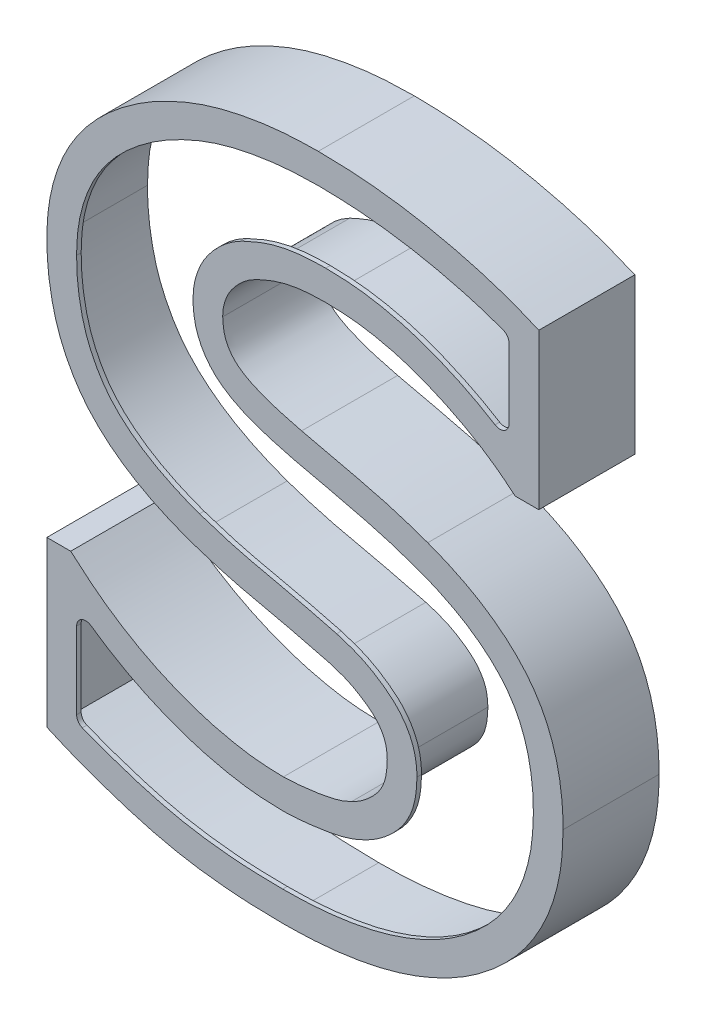
SolidWorks part; units mm, degrees
ref_plane "Front Plane" through (0, 0, 0) normal (0, 0, 1) x (1, 0, 0)
ref_plane "Top Plane" through (0, 0, 0) normal (0, 1, 0) x (1, 0, 0)
ref_plane "Right Plane" through (0, 0, 0) normal (1, 0, 0) x (0, 0, -1)
sketch "Sketch1" plane through (0, 0, 0) normal (0, 0, 1) x (1, 0, 0)
  line L30 (3196.1726, -1601.8231) -> (3190.9573, -1601.8231)
  line L31 (3190.9573, -1601.8231) -> (3190.9573, -1637.7551)
  line L32 (3293.3796, -1542.7978) -> (3298.5142, -1542.7978)
  line L33 (3298.5142, -1542.7978) -> (3298.5142, -1508.8154)
  line L34 (3196.1726, -1601.8231) -> (3190.9573, -1601.8231)
  line L35 (3190.9573, -1601.8231) -> (3190.9573, -1637.7551)
  line L36 (3293.3796, -1542.7978) -> (3298.5142, -1542.7978)
  line L37 (3298.5142, -1542.7978) -> (3298.5142, -1508.8154)
  spline S200 degree 3 poles (2284.4883, -3417.0637) (3101.6321, -1530.3936) (3137.0674, -1616.391) (3199.1425, -1641.1827) (3201.2322, -1641.9306) (3207.5334, -1644.0902) (3211.7766, -1645.3937) (3218.2649, -1646.912) (3220.4402, -1647.3415) (3224.8182, -1648.0349) (3227.02, -1648.3064) (3231.4398, -1648.7381) (3233.6526, -1648.8916) (3309.9762, -1651.9221) (3387.1158, -1589.7217) (3365.8768, -3641.246) knots -3.516933 -3.516933 -3.516933 -3.516933 0.125 0.125 0.25 0.25 0.5 0.5 0.625 0.625 0.75 0.75 0.875 0.875 5.055555 5.055555 5.055555 5.055555 only from (3190.9573, -1637.7551) to (3242.5214, -1649.127)
  spline S201 degree 3 poles (3389.1298, -3640.6843) (3110.4417, -1592.1851) (3184.4247, -1651.7096) (3249.8142, -1648.9185) (3251.6233, -1648.782) (3255.2229, -1648.3977) (3257.0144, -1648.156) (3260.5794, -1647.5655) (3262.3525, -1647.2137) (3265.8753, -1646.3706) (3267.6249, -1645.8785) (3270.2292, -1645.02) (3271.094, -1644.7142) (3272.8171, -1644.0635) (3273.6753, -1643.7187) (3277.9055, -1641.9116) (3281.1295, -1640.1881) (3284.9037, -1637.5903) (3285.6462, -1637.0493) (3287.1067, -1635.9249) (3287.8266, -1635.34) (3289.9254, -1633.5407) (3291.2507, -1632.2786) (3293.1156, -1630.2814) (3293.7161, -1629.5978) (3294.8692, -1628.1901) (3295.4216, -1627.4658) (3296.4798, -1625.9778) (3296.9856, -1625.2142) (3297.7103, -1624.0399) (3297.9462, -1623.6436) (3298.406, -1622.841) (3298.6305, -1622.4339) (3300.5824, -1618.7497) (3301.837, -1615.3159) (3302.8612, -1610.8435) (3303.0392, -1609.9402) (3303.3388, -1608.1148) (3303.46, -1607.1934) (3308.2244, -1558.5141) (3225.7698, -1504.7209) (5302.068, -1600.4559) knots -2.12183 -2.12183 -2.12183 -2.12183 0.0625 0.0625 0.125 0.125 0.1875 0.1875 0.25 0.25 0.3125 0.3125 0.34375 0.34375 0.375 0.375 0.5 0.5 0.53125 0.53125 0.5625 0.5625 0.625 0.625 0.65625 0.65625 0.6875 0.6875 0.71875 0.71875 0.734375 0.734375 0.75 0.75 0.875 0.875 0.90625 0.90625 0.9375 0.9375 2.557783 2.557783 2.557783 2.557783 only from (3242.5214, -1649.127) to (3303.831, -1600.7277)
  spline S202 degree 3 poles (5295.4273, -1434.3181) (3252.5035, -1691.2709) (3305.9059, -1640.2516) (3303.6811, -1596.2894) (3303.5852, -1595.1884) (3303.3185, -1592.9975) (3303.1491, -1591.9073) (3302.7301, -1589.7387) (3302.4809, -1588.6602) (3301.8832, -1586.5179) (3301.5302, -1585.4499) (3300.7417, -1583.3656) (3300.3092, -1582.3439) (3299.3308, -1580.3609) (3298.7826, -1579.4008) (3297.5897, -1577.5322) (3296.944, -1576.6227) (3295.5401, -1574.8697) (3294.7962, -1574.0388) (3293.2494, -1572.4406) (3292.4435, -1571.6767) (3290.7619, -1570.2245) (3289.8884, -1569.5338) (3288.0902, -1568.2079) (3287.165, -1567.5724) (3285.2879, -1566.3692) (3284.3308, -1565.8042) (3282.3786, -1564.749) (3281.3871, -1564.2518) (3279.3905, -1563.284) (3278.3817, -1562.8209) (3236.9653, -1545.6534) (3171.5196, -1578.3047) (4062.8736, 275.1184) knots -2.357405 -2.357405 -2.357405 -2.357405 0.0625 0.0625 0.125 0.125 0.1875 0.1875 0.25 0.25 0.3125 0.3125 0.375 0.375 0.4375 0.4375 0.5 0.5 0.5625 0.5625 0.625 0.625 0.6875 0.6875 0.75 0.75 0.8125 0.8125 0.875 0.875 0.9375 0.9375 3.393884 3.393884 3.393884 3.393884 only from (3303.831, -1600.7277) to (3274.2386, -1561.1811)
  spline S203 degree 3 poles (4092.8304, 259.838) (3375.1728, -1671.7225) (3333.4144, -1579.0951) (3265.1867, -1558.2212) (3262.8828, -1557.6217) (3129.3776, -1524.546) (2980.9575, -1565.3864) (3312.176, 431.8811) knots -6.989622 -6.989622 -6.989622 -6.989622 0.25 0.25 0.5 0.5 14.691826 14.691826 14.691826 14.691826 only from (3274.2386, -1561.1811) to (3246.6628, -1553.7945)
  spline S204 degree 3 poles (2866.7936, -3515.1405) (3367.7887, -1504.5868) (3293.2475, -1568.5546) (3240.5076, -1552.1032) (3240.0403, -1551.9495) (3239.115, -1551.6209) (3238.6566, -1551.4466) (3237.2855, -1550.9138) (3236.3715, -1550.5583) (3235.0513, -1549.905) (3234.6175, -1549.6684) (3233.7739, -1549.1585) (3233.3636, -1548.8885) (3232.5815, -1548.2976) (3232.2143, -1547.9707) (3231.5327, -1547.2476) (3231.2261, -1546.8629) (3230.6793, -1546.0529) (3230.4393, -1545.6268) (3230.1372, -1544.9511) (3230.0459, -1544.7184) (3229.8854, -1544.2495) (3229.8158, -1544.0128) (3229.6368, -1543.2965) (3229.5604, -1542.81) (3227.1802, -1519.9184) (3271.8943, -1489.2689) (1264.7707, -1913.0598) knots -6.715983 -6.715983 -6.715983 -6.715983 0.25 0.25 0.3125 0.3125 0.375 0.375 0.5 0.5 0.5625 0.5625 0.625 0.625 0.6875 0.6875 0.75 0.75 0.8125 0.8125 0.84375 0.84375 0.875 0.875 0.9375 0.9375 3.784326 3.784326 3.784326 3.784326 only from (3246.6628, -1553.7945) to (3229.4016, -1540.8359)
  spline S205 degree 3 poles (1256.17, -1216.6997) (3292.1305, -1587.2024) (3226.8255, -1556.6811) (3229.608, -1538.5806) (3229.7633, -1538.0366) (3230.1273, -1536.9587) (3230.3401, -1536.4237) (3230.8672, -1535.4276) (3231.1794, -1534.9602) (3231.8535, -1534.0569) (3232.219, -1533.6196) (3232.9898, -1532.7902) (3233.3942, -1532.3985) (3234.2421, -1531.6625) (3234.6849, -1531.3174) (3252.071, -1519.9003) (3307.7712, -1555.2808) (1935.0269, -12.1373) knots -3.809715 -3.809715 -3.809715 -3.809715 0.125 0.125 0.25 0.25 0.375 0.375 0.5 0.5 0.625 0.625 0.75 0.75 0.875 0.875 5.35521 5.35521 5.35521 5.35521 only from (3229.4016, -1540.8359) to (3236.6313, -1530.151)
  spline S206 degree 3 poles (2361.3876, 266.9714) (3202.1122, -1627.3675) (3205.7112, -1541.37) (3240.8796, -1528.3634) (3241.5073, -1528.1601) (3242.7729, -1527.8032) (3243.412, -1527.6489) (3244.7017, -1527.3856) (3245.3531, -1527.2765) (3246.6564, -1527.1014) (3247.3096, -1527.0353) (3288.8693, -1524.0388) (3334.8945, -1591.3649) (3225.703, 471.7079) knots -6.735966 -6.735966 -6.735966 -6.735966 0.25 0.25 0.375 0.375 0.5 0.5 0.625 0.625 0.75 0.75 8.561286 8.561286 8.561286 8.561286 only from (3236.6313, -1530.151) to (3251.9021, -1526.8487)
  spline S207 degree 3 poles (3313.4414, 470.4497) (3150.8906, -1604.2119) (3208.6341, -1522.6138) (3259.4657, -1527.2868) (3261.3369, -1527.5899) (3265.0638, -1528.346) (3266.9046, -1528.7955) (3270.5082, -1529.8837) (3272.2727, -1530.5241) (3275.7551, -1531.9257) (3277.4738, -1532.6845) (3280.0114, -1533.9274) (3280.8503, -1534.3596) (3282.5149, -1535.2582) (3283.3418, -1535.7253) (3285.7918, -1537.167) (3287.3889, -1538.1798) (3328.6344, -1568.0781) (3323.1117, -1661.3324) (4554.1151, 7.4638) knots -3.121892 -3.121892 -3.121892 -3.121892 0.125 0.125 0.25 0.25 0.375 0.375 0.5 0.5 0.625 0.625 0.6875 0.6875 0.75 0.75 0.875 0.875 4.120396 4.120396 4.120396 4.120396 only from (3251.9021, -1526.8487) to (3293.3796, -1542.7978)
  spline S208 degree 3 poles (4155.0848, 295.5208) (3380.8302, -1611.2773) (3348.4707, -1527.5834) (3290.8528, -1505.7529) (3288.8937, -1505.1035) (3284.9399, -1503.9045) (3282.9498, -1503.357) (3278.9444, -1502.3631) (3276.9288, -1501.9158) (3272.8794, -1501.1) (3270.8483, -1500.7338) (3266.7682, -1500.1188) (3264.7191, -1499.8687) (3260.6084, -1499.4578) (3258.5507, -1499.2984) (3189.0702, -1496.0526) (3118.2111, -1559.6931) (3156.4587, 495.3281) knots -3.48481 -3.48481 -3.48481 -3.48481 0.125 0.125 0.25 0.25 0.375 0.375 0.5 0.5 0.625 0.625 0.75 0.75 0.875 0.875 4.964131 4.964131 4.964131 4.964131 only from (3298.5142, -1508.8154) to (3250.3006, -1499.0381)
  spline S209 degree 3 poles (3057.6518, 488.9751) (3375.8631, -1556.8631) (3304.5949, -1496.2752) (3243.3298, -1499.2694) (3241.6033, -1499.4151) (3238.1713, -1499.8194) (3236.4652, -1500.0752) (3233.0727, -1500.693) (3231.386, -1501.0538) (3228.0358, -1501.9006) (3226.3729, -1502.3895) (3223.8996, -1503.2377) (3223.0787, -1503.5391) (3221.4439, -1504.1808) (3220.6281, -1504.5222) (3219.0159, -1505.2362) (3218.2192, -1505.6086) (3216.6427, -1506.381) (3215.8627, -1506.7806) (3214.3219, -1507.6115) (3213.5614, -1508.043) (3212.0631, -1508.9434) (3211.3258, -1509.413) (3209.8733, -1510.3881) (3209.158, -1510.8936) (3207.7477, -1511.9379) (3207.0524, -1512.4762) (3205.6844, -1513.5898) (3205.0106, -1514.1664) (3203.7034, -1515.3496) (3203.0687, -1515.9574) (3201.223, -1517.8307) (3200.0702, -1519.1462) (3198.4685, -1521.2285) (3197.9558, -1521.9409) (3197.2208, -1523.0385) (3196.9815, -1523.4093) (3196.5147, -1524.1609) (3196.287, -1524.5423) (3195.188, -1526.4602) (3194.4327, -1528.0404) (3193.1473, -1531.284) (3192.6145, -1532.9465) (3191.9738, -1535.499) (3191.7863, -1536.3595) (3191.4689, -1538.1017) (3191.3405, -1538.9764) (3186.4302, -1584.1219) (3271.7244, -1635.9395) (1192.8306, -1506.4458) knots -2.078551 -2.078551 -2.078551 -2.078551 0.0625 0.0625 0.125 0.125 0.1875 0.1875 0.25 0.25 0.3125 0.3125 0.34375 0.34375 0.375 0.375 0.40625 0.40625 0.4375 0.4375 0.46875 0.46875 0.5 0.5 0.53125 0.53125 0.5625 0.5625 0.59375 0.59375 0.625 0.625 0.6875 0.6875 0.71875 0.71875 0.734375 0.734375 0.75 0.75 0.8125 0.8125 0.875 0.875 0.90625 0.90625 0.9375 0.9375 2.51497 2.51497 2.51497 2.51497 only from (3250.3006, -1499.0381) to (3190.9569, -1545.139)
  spline S210 degree 3 poles (1201.1392, -1732.0358) (3244.5174, -1452.7478) (3188.7533, -1505.289) (3191.1209, -1549.8167) (3191.2265, -1550.9759) (3191.5206, -1553.2812) (3191.7095, -1554.4272) (3192.1555, -1556.7085) (3192.4102, -1557.8441) (3192.88, -1559.5337) (3193.0516, -1560.0945) (3193.4213, -1561.212) (3193.6197, -1561.7697) (3194.2435, -1563.4242) (3194.7001, -1564.5048) (3195.4775, -1566.0745) (3195.7509, -1566.59) (3196.3188, -1567.6091) (3196.6125, -1568.1133) (3197.2186, -1569.1113) (3197.5323, -1569.6045) (3198.191, -1570.5736) (3198.5371, -1571.0488) (3199.2623, -1571.9812) (3199.6411, -1572.439) (3200.415, -1573.3305) (3200.8108, -1573.7663) (3202.0258, -1575.0429) (3202.8738, -1575.8511) (3204.6443, -1577.384) (3205.5653, -1578.1103) (3207.467, -1579.4959) (3208.4501, -1580.1578) (3211.4486, -1582.033) (3213.5244, -1583.1254) (3216.7104, -1584.6157) (3217.786, -1585.0845) (3265.2111, -1604.2459) (3333.6583, -1577.5698) (2480.8499, -3442.3135) knots -2.261587 -2.261587 -2.261587 -2.261587 0.0625 0.0625 0.125 0.125 0.1875 0.1875 0.25 0.25 0.28125 0.28125 0.3125 0.3125 0.375 0.375 0.40625 0.40625 0.4375 0.4375 0.46875 0.46875 0.5 0.5 0.53125 0.53125 0.5625 0.5625 0.625 0.625 0.6875 0.6875 0.75 0.75 0.875 0.875 0.9375 0.9375 3.595499 3.595499 3.595499 3.595499 only from (3190.9569, -1545.139) to (3222.1685, -1586.7952)
  spline S211 degree 3 poles (2440.278, -3423.7139) (3120.3189, -1471.721) (3162.5464, -1570.4335) (3232.1823, -1589.8298) (3234.7307, -1590.4204) (3239.8366, -1591.564) (3242.3939, -1592.1176) (3331.9878, -1613.3076) (3404.2423, -1695.9129) (3964.6644, 267.953) knots -6.405604 -6.405604 -6.405604 -6.405604 0.25 0.25 0.5 0.5 0.75 0.75 9.298536 9.298536 9.298536 9.298536 only from (3222.1685, -1586.7952) to (3252.5513, -1594.6323)
  spline S212 degree 3 poles (3995.5228, 261.2808) (3149.9276, -1660.149) (3224.9032, -1581.6196) (3257.3722, -1596.3765) (3257.7242, -1596.5516) (3258.4164, -1596.9273) (3258.7572, -1597.1267) (3259.4319, -1597.5407) (3259.766, -1597.7545) (3260.4296, -1598.1925) (3260.7596, -1598.4186) (3261.7224, -1599.1248) (3262.3258, -1599.6356) (3263.1416, -1600.4949) (3263.3989, -1600.7964) (3263.8786, -1601.4359) (3264.1003, -1601.7737) (3264.4894, -1602.4677) (3264.6583, -1602.8265) (3264.9421, -1603.5693) (3265.0579, -1603.9562) (3265.2254, -1604.7412) (3265.2753, -1605.1376) (3267.1662, -1626.5474) (3227.8723, -1652.4053) (5257.5019, -1434.5975) knots -5.359923 -5.359923 -5.359923 -5.359923 0.25 0.25 0.3125 0.3125 0.375 0.375 0.4375 0.4375 0.5 0.5 0.625 0.625 0.6875 0.6875 0.75 0.75 0.8125 0.8125 0.875 0.875 0.9375 0.9375 4.235455 4.235455 4.235455 4.235455 only from (3252.5513, -1594.6323) to (3265.386, -1606.7339)
  spline S213 degree 3 poles (5253.2094, -1821.6114) (3168.1072, -1542.5744) (3271.3551, -1584.5463) (3264.9007, -1610.7395) (3264.8105, -1611.0404) (3264.5962, -1611.6351) (3264.4747, -1611.924) (3264.0743, -1612.7692) (3263.7625, -1613.306) (3263.0327, -1614.3163) (3262.604, -1614.7872) (3261.7186, -1615.6777) (3261.2626, -1616.1063) (3260.2999, -1616.9001) (3259.7919, -1617.2636) (3239.5943, -1629.7177) (3183.3286, -1596.203) (4528.1427, -3162.6322) knots -5.096482 -5.096482 -5.096482 -5.096482 0.25 0.25 0.3125 0.3125 0.375 0.375 0.5 0.5 0.625 0.625 0.75 0.75 0.875 0.875 5.469506 5.469506 5.469506 5.469506 only from (3265.386, -1606.7339) to (3257.5997, -1618.5148)
  spline S214 degree 3 poles (3885.0782, -3517.1586) (3277.2894, -1540.4289) (3276.0123, -1611.7526) (3255.2518, -1619.5179) (3254.6435, -1619.6966) (3253.4155, -1620.0156) (3252.795, -1620.1533) (3251.5459, -1620.4012) (3250.9164, -1620.5107) (3249.6536, -1620.7039) (3249.0206, -1620.7877) (3247.7527, -1620.9418) (3247.118, -1621.0135) (3245.8471, -1621.142) (3245.2113, -1621.2001) (3214.9983, -1623.1368) (3182.2112, -1575.7571) (3285.7343, -3620.1449) knots -4.109234 -4.109234 -4.109234 -4.109234 0.125 0.125 0.25 0.25 0.375 0.375 0.5 0.5 0.625 0.625 0.75 0.75 0.875 0.875 6.679038 6.679038 6.679038 6.679038 only from (3257.5997, -1618.5148) to (3242.6603, -1621.3162)
  spline S215 degree 3 poles (3142.4723, -3617.0203) (3341.9672, -1578.2296) (3287.7888, -1623.6098) (3238.3507, -1621.1495) (3237.2778, -1621.071) (3235.143, -1620.8233) (3234.0805, -1620.6591) (3231.9624, -1620.2746) (3230.9066, -1620.0557) (3228.7998, -1619.578) (3227.7515, -1619.3172) (3225.6786, -1618.7481) (3224.6527, -1618.4385) (3221.6069, -1617.4342) (3219.6167, -1616.6691) (3215.7004, -1614.9871) (3213.7767, -1614.0645) (3210.9494, -1612.5428) (3210.0163, -1612.0133) (3208.1677, -1610.9128) (3207.2505, -1610.3411) (3204.5409, -1608.5756) (3202.7905, -1607.3254) (3154.4905, -1568.8851) (3152.7107, -1473.2001) (1849.9523, -3077.3406) knots -2.746767 -2.746767 -2.746767 -2.746767 0.0625 0.0625 0.125 0.125 0.1875 0.1875 0.25 0.25 0.3125 0.3125 0.375 0.375 0.5 0.5 0.625 0.625 0.6875 0.6875 0.75 0.75 0.875 0.875 4.338516 4.338516 4.338516 4.338516 only from (3242.6603, -1621.3162) to (3196.1726, -1601.8231)
  spline S216 degree 3 poles (3190.9573, -1637.7551) (3192.9918, -1638.6416) (3195.0227, -1639.5373) (3199.1425, -1641.1827) (3201.2322, -1641.9306) (3207.5334, -1644.0902) (3211.7766, -1645.3937) (3218.2649, -1646.912) (3220.4402, -1647.3415) (3224.8182, -1648.0349) (3227.02, -1648.3064) (3231.4398, -1648.7381) (3233.6526, -1648.8916) (3238.0843, -1649.0675) (3240.3029, -1649.0973) (3242.5214, -1649.127) knots 0 0 0 0 0.125 0.125 0.25 0.25 0.5 0.5 0.625 0.625 0.75 0.75 0.875 0.875 1 1 1 1
  spline S217 degree 3 poles (3242.5214, -1649.127) (3244.3489, -1649.1005) (3246.1764, -1649.0738) (3249.8142, -1648.9185) (3251.6233, -1648.782) (3255.2229, -1648.3977) (3257.0144, -1648.156) (3260.5794, -1647.5655) (3262.3525, -1647.2137) (3265.8753, -1646.3706) (3267.6249, -1645.8785) (3270.2292, -1645.02) (3271.094, -1644.7142) (3272.8171, -1644.0635) (3273.6753, -1643.7187) (3277.9055, -1641.9116) (3281.1295, -1640.1881) (3284.9037, -1637.5903) (3285.6462, -1637.0493) (3287.1067, -1635.9249) (3287.8266, -1635.34) (3289.9254, -1633.5407) (3291.2507, -1632.2786) (3293.1156, -1630.2814) (3293.7161, -1629.5978) (3294.8692, -1628.1901) (3295.4216, -1627.4658) (3296.4798, -1625.9778) (3296.9856, -1625.2142) (3297.7103, -1624.0399) (3297.9462, -1623.6436) (3298.406, -1622.841) (3298.6305, -1622.4339) (3300.5824, -1618.7497) (3301.837, -1615.3159) (3302.8612, -1610.8435) (3303.0392, -1609.9402) (3303.3388, -1608.1148) (3303.46, -1607.1934) (3303.7305, -1604.4301) (3303.7811, -1602.5789) (3303.831, -1600.7277) knots 0 0 0 0 0.0625 0.0625 0.125 0.125 0.1875 0.1875 0.25 0.25 0.3125 0.3125 0.34375 0.34375 0.375 0.375 0.5 0.5 0.53125 0.53125 0.5625 0.5625 0.625 0.625 0.65625 0.65625 0.6875 0.6875 0.71875 0.71875 0.734375 0.734375 0.75 0.75 0.875 0.875 0.90625 0.90625 0.9375 0.9375 1 1 1 1
  spline S218 degree 3 poles (3303.831, -1600.7277) (3303.8121, -1599.6154) (3303.7931, -1598.5031) (3303.6811, -1596.2894) (3303.5852, -1595.1884) (3303.3185, -1592.9975) (3303.1491, -1591.9073) (3302.7301, -1589.7387) (3302.4809, -1588.6602) (3301.8832, -1586.5179) (3301.5302, -1585.4499) (3300.7417, -1583.3656) (3300.3092, -1582.3439) (3299.3308, -1580.3609) (3298.7826, -1579.4008) (3297.5897, -1577.5322) (3296.944, -1576.6227) (3295.5401, -1574.8697) (3294.7962, -1574.0388) (3293.2494, -1572.4406) (3292.4435, -1571.6767) (3290.7619, -1570.2245) (3289.8884, -1569.5338) (3288.0902, -1568.2079) (3287.165, -1567.5724) (3285.2879, -1566.3692) (3284.3308, -1565.8042) (3282.3786, -1564.749) (3281.3871, -1564.2518) (3279.3905, -1563.284) (3278.3817, -1562.8209) (3276.3264, -1561.969) (3275.2825, -1561.575) (3274.2386, -1561.1811) knots 0 0 0 0 0.0625 0.0625 0.125 0.125 0.1875 0.1875 0.25 0.25 0.3125 0.3125 0.375 0.375 0.4375 0.4375 0.5 0.5 0.5625 0.5625 0.625 0.625 0.6875 0.6875 0.75 0.75 0.8125 0.8125 0.875 0.875 0.9375 0.9375 1 1 1 1
  spline S219 degree 3 poles (3274.2386, -1561.1811) (3271.9901, -1560.3979) (3269.7415, -1559.6147) (3265.1867, -1558.2212) (3262.8828, -1557.6217) (3255.9496, -1555.904) (3251.306, -1554.8499) (3246.6628, -1553.7945) knots 0 0 0 0 0.25 0.25 0.5 0.5 1 1 1 1
  spline S220 degree 3 poles (3246.6628, -1553.7945) (3244.7572, -1553.3165) (3242.8525, -1552.8347) (3240.5076, -1552.1032) (3240.0403, -1551.9495) (3239.115, -1551.6209) (3238.6566, -1551.4466) (3237.2855, -1550.9138) (3236.3715, -1550.5583) (3235.0513, -1549.905) (3234.6175, -1549.6684) (3233.7739, -1549.1585) (3233.3636, -1548.8885) (3232.5815, -1548.2976) (3232.2143, -1547.9707) (3231.5327, -1547.2476) (3231.2261, -1546.8629) (3230.6793, -1546.0529) (3230.4393, -1545.6268) (3230.1372, -1544.9511) (3230.0459, -1544.7184) (3229.8854, -1544.2495) (3229.8158, -1544.0128) (3229.6368, -1543.2965) (3229.5604, -1542.81) (3229.4581, -1541.8265) (3229.4296, -1541.3307) (3229.4016, -1540.8359) knots 0 0 0 0 0.25 0.25 0.3125 0.3125 0.375 0.375 0.5 0.5 0.5625 0.5625 0.625 0.625 0.6875 0.6875 0.75 0.75 0.8125 0.8125 0.84375 0.84375 0.875 0.875 0.9375 0.9375 1 1 1 1
  spline S221 degree 3 poles (3229.4016, -1540.8359) (3229.4196, -1540.2657) (3229.4367, -1539.6953) (3229.608, -1538.5806) (3229.7633, -1538.0366) (3230.1273, -1536.9587) (3230.3401, -1536.4237) (3230.8672, -1535.4276) (3231.1794, -1534.9602) (3231.8535, -1534.0569) (3232.219, -1533.6196) (3232.9898, -1532.7902) (3233.3942, -1532.3985) (3234.2421, -1531.6625) (3234.6849, -1531.3174) (3235.6288, -1530.6976) (3236.1309, -1530.4239) (3236.6313, -1530.151) knots 0 0 0 0 0.125 0.125 0.25 0.25 0.375 0.375 0.5 0.5 0.625 0.625 0.75 0.75 0.875 0.875 1 1 1 1
  spline S222 degree 3 poles (3236.6313, -1530.151) (3237.8282, -1529.6003) (3239.025, -1529.0493) (3240.8796, -1528.3634) (3241.5073, -1528.1601) (3242.7729, -1527.8032) (3243.412, -1527.6489) (3244.7017, -1527.3856) (3245.3531, -1527.2765) (3246.6564, -1527.1014) (3247.3096, -1527.0353) (3249.2733, -1526.8937) (3250.5877, -1526.8713) (3251.9021, -1526.8487) knots 0 0 0 0 0.25 0.25 0.375 0.375 0.5 0.5 0.625 0.625 0.75 0.75 1 1 1 1
  spline S223 degree 3 poles (3251.9021, -1526.8487) (3253.7995, -1526.8947) (3255.697, -1526.9403) (3259.4657, -1527.2868) (3261.3369, -1527.5899) (3265.0638, -1528.346) (3266.9046, -1528.7955) (3270.5082, -1529.8837) (3272.2727, -1530.5241) (3275.7551, -1531.9257) (3277.4738, -1532.6845) (3280.0114, -1533.9274) (3280.8503, -1534.3596) (3282.5149, -1535.2582) (3283.3418, -1535.7253) (3285.7918, -1537.167) (3287.3889, -1538.1798) (3290.4483, -1540.3975) (3291.9109, -1541.602) (3293.3796, -1542.7978) knots 0 0 0 0 0.125 0.125 0.25 0.25 0.375 0.375 0.5 0.5 0.625 0.625 0.6875 0.6875 0.75 0.75 0.875 0.875 1 1 1 1
  spline S224 degree 3 poles (3298.5142, -1508.8154) (3296.61, -1508.0199) (3294.7096, -1507.2142) (3290.8528, -1505.7529) (3288.8937, -1505.1035) (3284.9399, -1503.9045) (3282.9498, -1503.357) (3278.9444, -1502.3631) (3276.9288, -1501.9158) (3272.8794, -1501.1) (3270.8483, -1500.7338) (3266.7682, -1500.1188) (3264.7191, -1499.8687) (3260.6084, -1499.4578) (3258.5507, -1499.2984) (3254.4289, -1499.1058) (3252.3647, -1499.0719) (3250.3006, -1499.0381) knots 0 0 0 0 0.125 0.125 0.25 0.25 0.375 0.375 0.5 0.5 0.625 0.625 0.75 0.75 0.875 0.875 1 1 1 1
  spline S225 degree 3 poles (3250.3006, -1499.0381) (3248.5529, -1499.0687) (3246.8052, -1499.0996) (3243.3298, -1499.2694) (3241.6033, -1499.4151) (3238.1713, -1499.8194) (3236.4652, -1500.0752) (3233.0727, -1500.693) (3231.386, -1501.0538) (3228.0358, -1501.9006) (3226.3729, -1502.3895) (3223.8996, -1503.2377) (3223.0787, -1503.5391) (3221.4439, -1504.1808) (3220.6281, -1504.5222) (3219.0159, -1505.2362) (3218.2192, -1505.6086) (3216.6427, -1506.381) (3215.8627, -1506.7806) (3214.3219, -1507.6115) (3213.5614, -1508.043) (3212.0631, -1508.9434) (3211.3258, -1509.413) (3209.8733, -1510.3881) (3209.158, -1510.8936) (3207.7477, -1511.9379) (3207.0524, -1512.4762) (3205.6844, -1513.5898) (3205.0106, -1514.1664) (3203.7034, -1515.3496) (3203.0687, -1515.9574) (3201.223, -1517.8307) (3200.0702, -1519.1462) (3198.4685, -1521.2285) (3197.9558, -1521.9409) (3197.2208, -1523.0385) (3196.9815, -1523.4093) (3196.5147, -1524.1609) (3196.287, -1524.5423) (3195.188, -1526.4602) (3194.4327, -1528.0404) (3193.1473, -1531.284) (3192.6145, -1532.9465) (3191.9738, -1535.499) (3191.7863, -1536.3595) (3191.4689, -1538.1017) (3191.3405, -1538.9764) (3191.0543, -1541.6073) (3191.005, -1543.3731) (3190.9569, -1545.139) knots 0 0 0 0 0.0625 0.0625 0.125 0.125 0.1875 0.1875 0.25 0.25 0.3125 0.3125 0.34375 0.34375 0.375 0.375 0.40625 0.40625 0.4375 0.4375 0.46875 0.46875 0.5 0.5 0.53125 0.53125 0.5625 0.5625 0.59375 0.59375 0.625 0.625 0.6875 0.6875 0.71875 0.71875 0.734375 0.734375 0.75 0.75 0.8125 0.8125 0.875 0.875 0.90625 0.90625 0.9375 0.9375 1 1 1 1
  spline S226 degree 3 poles (3190.9569, -1545.139) (3190.9769, -1546.3118) (3190.9969, -1547.4845) (3191.1209, -1549.8167) (3191.2265, -1550.9759) (3191.5206, -1553.2812) (3191.7095, -1554.4272) (3192.1555, -1556.7085) (3192.4102, -1557.8441) (3192.88, -1559.5337) (3193.0516, -1560.0945) (3193.4213, -1561.212) (3193.6197, -1561.7697) (3194.2435, -1563.4242) (3194.7001, -1564.5048) (3195.4775, -1566.0745) (3195.7509, -1566.59) (3196.3188, -1567.6091) (3196.6125, -1568.1133) (3197.2186, -1569.1113) (3197.5323, -1569.6045) (3198.191, -1570.5736) (3198.5371, -1571.0488) (3199.2623, -1571.9812) (3199.6411, -1572.439) (3200.415, -1573.3305) (3200.8108, -1573.7663) (3202.0258, -1575.0429) (3202.8738, -1575.8511) (3204.6443, -1577.384) (3205.5653, -1578.1103) (3207.467, -1579.4959) (3208.4501, -1580.1578) (3211.4486, -1582.033) (3213.5244, -1583.1254) (3216.7104, -1584.6157) (3217.786, -1585.0845) (3219.9651, -1585.9649) (3221.0668, -1586.38) (3222.1685, -1586.7952) knots 0 0 0 0 0.0625 0.0625 0.125 0.125 0.1875 0.1875 0.25 0.25 0.28125 0.28125 0.3125 0.3125 0.375 0.375 0.40625 0.40625 0.4375 0.4375 0.46875 0.46875 0.5 0.5 0.53125 0.53125 0.5625 0.5625 0.625 0.625 0.6875 0.6875 0.75 0.75 0.875 0.875 0.9375 0.9375 1 1 1 1
  spline S227 degree 3 poles (3222.1685, -1586.7952) (3224.6544, -1587.6103) (3227.1403, -1588.4254) (3232.1823, -1589.8298) (3234.7307, -1590.4204) (3239.8366, -1591.564) (3242.3939, -1592.1176) (3247.4853, -1593.3218) (3250.0183, -1593.9769) (3252.5513, -1594.6323) knots 0 0 0 0 0.25 0.25 0.5 0.5 0.75 0.75 1 1 1 1
  spline S228 degree 3 poles (3252.5513, -1594.6323) (3254.0673, -1595.0981) (3255.5834, -1595.5635) (3257.3722, -1596.3765) (3257.7242, -1596.5516) (3258.4164, -1596.9273) (3258.7572, -1597.1267) (3259.4319, -1597.5407) (3259.766, -1597.7545) (3260.4296, -1598.1925) (3260.7596, -1598.4186) (3261.7224, -1599.1248) (3262.3258, -1599.6356) (3263.1416, -1600.4949) (3263.3989, -1600.7964) (3263.8786, -1601.4359) (3264.1003, -1601.7737) (3264.4894, -1602.4677) (3264.6583, -1602.8265) (3264.9421, -1603.5693) (3265.0579, -1603.9562) (3265.2254, -1604.7412) (3265.2753, -1605.1376) (3265.3457, -1605.934) (3265.3661, -1606.334) (3265.386, -1606.7339) knots 0 0 0 0 0.25 0.25 0.3125 0.3125 0.375 0.375 0.4375 0.4375 0.5 0.5 0.625 0.625 0.6875 0.6875 0.75 0.75 0.8125 0.8125 0.875 0.875 0.9375 0.9375 1 1 1 1
  spline S229 degree 3 poles (3265.386, -1606.7339) (3265.3322, -1607.9804) (3265.2736, -1609.2262) (3264.9007, -1610.7395) (3264.8105, -1611.0404) (3264.5962, -1611.6351) (3264.4747, -1611.924) (3264.0743, -1612.7692) (3263.7625, -1613.306) (3263.0327, -1614.3163) (3262.604, -1614.7872) (3261.7186, -1615.6777) (3261.2626, -1616.1063) (3260.2999, -1616.9001) (3259.7919, -1617.2636) (3258.722, -1617.9233) (3258.1599, -1618.2194) (3257.5997, -1618.5148) knots 0 0 0 0 0.25 0.25 0.3125 0.3125 0.375 0.375 0.5 0.5 0.625 0.625 0.75 0.75 0.875 0.875 1 1 1 1
  spline S230 degree 3 poles (3257.5997, -1618.5148) (3257.0213, -1618.7943) (3256.4424, -1619.0726) (3255.2518, -1619.5179) (3254.6435, -1619.6966) (3253.4155, -1620.0156) (3252.795, -1620.1533) (3251.5459, -1620.4012) (3250.9164, -1620.5107) (3249.6536, -1620.7039) (3249.0206, -1620.7877) (3247.7527, -1620.9418) (3247.118, -1621.0135) (3245.8471, -1621.142) (3245.2113, -1621.2001) (3243.9373, -1621.2817) (3243.2988, -1621.2997) (3242.6603, -1621.3162) knots 0 0 0 0 0.125 0.125 0.25 0.25 0.375 0.375 0.5 0.5 0.625 0.625 0.75 0.75 0.875 0.875 1 1 1 1
  spline S231 degree 3 poles (3242.6603, -1621.3162) (3241.5814, -1621.2865) (3240.5026, -1621.2566) (3238.3507, -1621.1495) (3237.2778, -1621.071) (3235.143, -1620.8233) (3234.0805, -1620.6591) (3231.9624, -1620.2746) (3230.9066, -1620.0557) (3228.7998, -1619.578) (3227.7515, -1619.3172) (3225.6786, -1618.7481) (3224.6527, -1618.4385) (3221.6069, -1617.4342) (3219.6167, -1616.6691) (3215.7004, -1614.9871) (3213.7767, -1614.0645) (3210.9494, -1612.5428) (3210.0163, -1612.0133) (3208.1677, -1610.9128) (3207.2505, -1610.3411) (3204.5409, -1608.5756) (3202.7905, -1607.3254) (3199.4256, -1604.6473) (3197.8016, -1603.232) (3196.1726, -1601.8231) knots 0 0 0 0 0.0625 0.0625 0.125 0.125 0.1875 0.1875 0.25 0.25 0.3125 0.3125 0.375 0.375 0.5 0.5 0.625 0.625 0.6875 0.6875 0.75 0.75 0.875 0.875 1 1 1 1
  dimension "D1" = 1.5
extrude "Boss-Extrude1" add sketch "Sketch1" along normal blind 1 and the other way blind 20
sketch3d "3DSketch3"
  line L0 (3197.4573, -1611.3857, 1) -> (3197.4573, -1633.4798, 1)
  line L1 (3292.0142, -1533.5232, 1) -> (3292.0142, -1513.1649, 1)
  line L2 (3197.4573, -1611.3857, 1) -> (3197.4573, -1633.4798, 1)
  line L3 (3292.0142, -1533.5232, 1) -> (3292.0142, -1513.1649, 1)
  spline S0 degree 5 poles (4580.7215, -263.8915, 1) (3283.2461, -1350.3751, 1) (3280.2183, -1414.0576, 1) (3277.4391, -1478.3768, 1) (3274.6532, -1542.8424, 1) (3271.8673, -1607.3079, 1) (3271.8608, -1607.4546, 1) (3271.8382, -1607.9355, 1) (3271.8097, -1608.4161, 1) (3271.786, -1608.7499, 1) (3271.7169, -1609.5582, 1) (3271.6132, -1610.3639, 1) (3271.5385, -1610.8353, 1) (3271.3594, -1611.7637, 1) (3271.1114, -1612.6761, 1) (3270.9719, -1613.1235, 1) (3270.6776, -1613.958, 1) (3270.3261, -1614.7697, 1) (3270.1487, -1615.1464, 1) (3269.7472, -1615.9347, 1) (3269.2967, -1616.6965, 1) (3269.0442, -1617.0909, 1) (3268.4933, -1617.8843, 1) (3267.8795, -1618.6301, 1) (3267.5495, -1619.0034, 1) (3266.8353, -1619.7667, 1) (3266.0881, -1620.4958, 1) (3265.6873, -1620.8665, 1) (3264.8931, -1621.5588, 1) (3264.056, -1622.2006, 1) (3263.6431, -1622.4975, 1) (3262.9387, -1622.9708, 1) (3262.2104, -1623.4047, 1) (3261.9153, -1623.5734, 1) (3261.4816, -1623.8132, 1) (3261.0445, -1624.0464, 1) (3260.9071, -1624.1191, 1) (3241.3524, -1634.4319, 1) (3221.7978, -1644.7447, 1) (3202.3811, -1654.9849, 1) (3181.9636, -1665.1517, 1) (5168.8746, -2021.4633, 1) knots -14.491372 -14.491372 -14.491372 -14.491372 -14.491372 -14.491372 0.013641 0.013641 0.013641 0.046719 0.046719 0.046719 0.122101 0.122101 0.122101 0.229433 0.229433 0.229433 0.334825 0.334825 0.334825 0.428531 0.428531 0.428531 0.533896 0.533896 0.533896 0.645937 0.645937 0.645937 0.768868 0.768868 0.768868 0.883239 0.883239 0.883239 0.959797 0.959797 0.959797 0.994843 0.994843 0.994843 5.940746 5.940746 5.940746 5.940746 5.940746 5.940746 only from (3271.8931, -1606.7121, 1) to (3260.5307, -1624.3177, 1)
  spline S1 degree 5 poles (3223.8625, -197.3996, 1.1184) (3343.4985, -1584.7595, 0.9999) (3322.9394, -1594.1627, 1) (3302.1021, -1604.2311, 1) (3281.0632, -1614.3967, 1) (3260.0242, -1624.5623, 1) (3259.8221, -1624.6589, 1) (3259.2208, -1624.94, 1) (3258.6083, -1625.1983, 1) (3258.1981, -1625.3592, 1) (3257.183, -1625.728, 1) (3256.148, -1626.0322, 1) (3255.5298, -1626.1937, 1) (3254.3212, -1626.4788, 1) (3253.1043, -1626.723, 1) (3252.512, -1626.8322, 1) (3251.3507, -1627.0282, 1) (3250.1845, -1627.1914, 1) (3249.6138, -1627.265, 1) (3248.481, -1627.4019, 1) (3247.347, -1627.5274, 1) (3246.7845, -1627.5851, 1) (3245.8453, -1627.6706, 1) (3244.904, -1627.7336, 1) (3244.5268, -1627.755, 1) (3243.9608, -1627.7815, 1) (3243.3945, -1627.7991, 1) (3243.2058, -1627.8043, 1) (3204.6966, -1628.7998, 1) (3166.1875, -1629.7953, 1) (3127.867, -1630.7861, 1) (3089.0792, -1631.1931, 1) (4934.0875, -2275.4629, 1) knots -6.300977 -6.300977 -6.300977 -6.300977 -6.300977 -6.300977 0.006238 0.006238 0.006238 0.067287 0.067287 0.067287 0.187111 0.187111 0.187111 0.361112 0.361112 0.361112 0.525229 0.525229 0.525229 0.682047 0.682047 0.682047 0.836146 0.836146 0.836146 0.939081 0.939081 0.939081 0.990541 0.990541 0.990541 11.437972 11.437972 11.437972 11.437972 11.437972 11.437972 only from (3260.5307, -1624.3177, 1) to (3242.6548, -1627.8185, 1)
  spline S2 degree 5 poles (4319.6493, -222.7025, 0.7374) (3399.7098, -1632.6519, 1.0002) (3360.7613, -1631.0716, 1) (3321.3345, -1629.9857, 1) (3281.5329, -1628.8894, 1) (3241.7314, -1627.7931, 1) (3241.3564, -1627.7823, 1) (3240.2368, -1627.7477, 1) (3239.1172, -1627.7016, 1) (3238.373, -1627.6627, 1) (3236.4973, -1627.5353, 1) (3234.6298, -1627.314, 1) (3233.5059, -1627.1506, 1) (3231.2673, -1626.7737, 1) (3229.0456, -1626.3142, 1) (3227.9403, -1626.0641, 1) (3225.7358, -1625.5222, 1) (3223.5525, -1624.8986, 1) (3222.465, -1624.5657, 1) (3220.1798, -1623.8181, 1) (3217.9274, -1622.9773, 1) (3216.7495, -1622.5098, 1) (3214.271, -1621.4695, 1) (3211.8351, -1620.3324, 1) (3210.5608, -1619.7039, 1) (3208.2246, -1618.4865, 1) (3205.942, -1617.1709, 1) (3204.902, -1616.5449, 1) (3203.1474, -1615.4449, 1) (3201.4273, -1614.2931, 1) (3200.7217, -1613.807, 1) (3153.3295, -1580.1787, 1) (3139.8774, -1499.8277, 1) (3313.3196, -1324.604, 1) (3827.2077, -1002.6208, 1) (4835.2681, -483.1895, 1) knots -4.027061 -4.027061 -4.027061 -4.027061 -4.027061 -4.027061 0.003547 0.003547 0.003547 0.04188 0.04188 0.04188 0.118001 0.118001 0.118001 0.233967 0.233967 0.233967 0.349743 0.349743 0.349743 0.465899 0.465899 0.465899 0.59535 0.59535 0.59535 0.740447 0.740447 0.740447 0.8644 0.8644 0.8644 0.951944 0.951944 0.951944 6.802332 6.802332 6.802332 6.802332 6.802332 6.802332 only from (3242.6548, -1627.8185, 1) to (3197.4573, -1611.3857, 1)
  spline S3 degree 5 poles (2341.4314, -3437.2251, 1) (2797.6514, -2285.0387, 1) (3036.5338, -1736.9031, 1) (3133.1938, -1584.6028, 1) (3163.8213, -1621.2041, 1) (3203.0537, -1635.6893, 1) (3204.4352, -1636.1744, 1) (3207.1943, -1637.1059, 1) (3209.9677, -1637.9919, 1) (3211.3511, -1638.4168, 1) (3214.104, -1639.2194, 1) (3216.8841, -1639.9275, 1) (3218.2677, -1640.2524, 1) (3221.0483, -1640.846, 1) (3223.852, -1641.316, 1) (3225.2592, -1641.5232, 1) (3228.1021, -1641.8906, 1) (3230.9547, -1642.1691, 1) (3232.3937, -1642.2861, 1) (3234.8079, -1642.442, 1) (3237.2252, -1642.5286, 1) (3238.2004, -1642.5549, 1) (3282.5446, -1643.4713, 1) (3326.8658, -1637.1017, 1) (3370.8401, -1828.8727, 1) (3416.0924, -2423.6137, 1) (3463.2695, -3626.2955, 1) knots -4.289829 -4.289829 -4.289829 -4.289829 -4.289829 -4.289829 0.066713 0.066713 0.066713 0.22474 0.22474 0.22474 0.38096 0.38096 0.38096 0.534292 0.534292 0.534292 0.687778 0.687778 0.687778 0.843593 0.843593 0.843593 0.948894 0.948894 0.948894 5.631235 5.631235 5.631235 5.631235 5.631235 5.631235 only from (3197.4573, -1633.4798, 1) to (3242.5177, -1642.6264, 1)
  spline S4 degree 5 poles (3045.4395, -3629.6288, 1) (3086.9335, -2427.6447, 1) (3127.1311, -1831.867, 1) (3166.4393, -1638.3815, 1) (3205.9968, -1643.353, 1) (3245.5671, -1642.5752, 1) (3246.255, -1642.5581, 1) (3247.9669, -1642.5021, 1) (3249.6771, -1642.4013, 1) (3250.6993, -1642.3251, 1) (3252.719, -1642.1434, 1) (3254.7323, -1641.9011, 1) (3255.7261, -1641.7665, 1) (3257.8106, -1641.4523, 1) (3259.8846, -1641.0725, 1) (3260.968, -1640.8531, 1) (3263.2302, -1640.3455, 1) (3265.4663, -1639.7283, 1) (3266.628, -1639.3755, 1) (3269.0186, -1638.5821, 1) (3271.3631, -1637.6615, 1) (3272.5634, -1637.1495, 1) (3274.8271, -1636.1022, 1) (3277.0251, -1634.9201, 1) (3278.0558, -1634.3246, 1) (3279.9689, -1633.1349, 1) (3281.7996, -1631.8235, 1) (3282.6449, -1631.1792, 1) (3284.2081, -1629.915, 1) (3285.7028, -1628.5704, 1) (3286.39, -1627.9179, 1) (3287.7175, -1626.5816, 1) (3288.9597, -1625.1643, 1) (3289.5542, -1624.4403, 1) (3290.6873, -1622.9625, 1) (3291.7163, -1621.4105, 1) (3292.2017, -1620.6222, 1) (3293.1231, -1619.0093, 1) (3293.9379, -1617.3401, 1) (3294.3189, -1616.4896, 1) (3294.9853, -1614.8578, 1) (3295.5456, -1613.1869, 1) (3295.7867, -1612.3916, 1) (3296.1978, -1610.8858, 1) (3296.5322, -1609.3618, 1) (3296.6711, -1608.6455, 1) (3296.8998, -1607.2811, 1) (3297.0597, -1605.9071, 1) (3297.1214, -1605.2559, 1) (3297.2039, -1604.1617, 1) (3297.2555, -1603.0661, 1) (3297.2725, -1602.6233, 1) (3298.2184, -1573.7513, 1) (3293.8964, -1544.7793, 1) (3488.7696, -1520.0305, 1) (4087.0085, -1502.9358, 1) (5292.8699, -1497.4605, 1) knots -2.483516 -2.483516 -2.483516 -2.483516 -2.483516 -2.483516 0.021561 0.021561 0.021561 0.06589 0.06589 0.06589 0.131897 0.131897 0.131897 0.196489 0.196489 0.196489 0.267667 0.267667 0.267667 0.3458 0.3458 0.3458 0.429771 0.429771 0.429771 0.506327 0.506327 0.506327 0.574732 0.574732 0.574732 0.635718 0.635718 0.635718 0.695982 0.695982 0.695982 0.755532 0.755532 0.755532 0.81548 0.81548 0.81548 0.868947 0.868947 0.868947 0.915915 0.915915 0.915915 0.958025 0.958025 0.958025 0.986568 0.986568 0.986568 2.818876 2.818876 2.818876 2.818876 2.818876 2.818876 only from (3242.5177, -1642.6264, 1) to (3297.3295, -1600.6954, 1)
  spline S5 degree 5 poles (5291.4165, -1733.4676, 1) (4086.2891, -1705.2371, 1) (3488.2595, -1678.1028, 1) (3293.462, -1651.7484, 1) (3297.901, -1625.3811, 1) (3297.2961, -1599.0041, 1) (3297.2847, -1598.6061, 1) (3297.2474, -1597.62, 1) (3297.1808, -1596.6352, 1) (3297.1307, -1596.0485, 1) (3297.012, -1594.8984, 1) (3296.8535, -1593.7533, 1) (3296.766, -1593.1927, 1) (3296.5725, -1592.0807, 1) (3296.3398, -1590.9759, 1) (3296.2132, -1590.4288, 1) (3295.9391, -1589.3509, 1) (3295.6141, -1588.2873, 1) (3295.4415, -1587.7641, 1) (3295.0787, -1586.7371, 1) (3294.6764, -1585.7246, 1) (3294.4662, -1585.229, 1) (3294.023, -1584.257, 1) (3293.5218, -1583.3132, 1) (3293.2597, -1582.8519, 1) (3292.6145, -1581.7849, 1) (3291.9061, -1580.7591, 1) (3291.4789, -1580.184, 1) (3290.4543, -1578.8987, 1) (3289.3316, -1577.6958, 1) (3288.6708, -1577.0424, 1) (3287.2926, -1575.7758, 1) (3285.8352, -1574.6055, 1) (3285.0832, -1574.0396, 1) (3283.6802, -1573.0466, 1) (3282.2304, -1572.1248, 1) (3281.565, -1571.7226, 1) (3280.3794, -1571.0422, 1) (3279.1678, -1570.4102, 1) (3278.6413, -1570.1449, 1) (3277.5653, -1569.6175, 1) (3276.4812, -1569.1068, 1) (3275.9277, -1568.8539, 1) (3274.9988, -1568.4467, 1) (3274.0575, -1568.0693, 1) (3273.6794, -1567.9218, 1) (3247.859, -1558.0255, 1) (3220.5104, -1552.705, 1) (3256.5455, -1358.8784, 1) (3420.0288, -783.4411, 1) (3775.3572, 366.5971, 1) knots -2.84576 -2.84576 -2.84576 -2.84576 -2.84576 -2.84576 0.019748 0.019748 0.019748 0.063657 0.063657 0.063657 0.128567 0.128567 0.128567 0.191118 0.191118 0.191118 0.253005 0.253005 0.253005 0.313731 0.313731 0.313731 0.373049 0.373049 0.373049 0.431494 0.431494 0.431494 0.510413 0.510413 0.510413 0.612582 0.612582 0.612582 0.716237 0.716237 0.716237 0.801931 0.801931 0.801931 0.866942 0.866942 0.866942 0.934043 0.934043 0.934043 0.97879 0.97879 0.97879 3.983026 3.983026 3.983026 3.983026 3.983026 3.983026 only from (3297.3295, -1600.6954, 1) to (3272.0218, -1567.292, 1)
  spline S6 degree 5 poles (4164.4802, 218.1482, 1) (3705.2809, -890.8014, 1) (3457.25, -1433.2692, 1) (3349.4466, -1599.7345, 1) (3310.169, -1580.3872, 1) (3268.9557, -1566.2304, 1) (3268.2706, -1565.9986, 1) (3266.5518, -1565.4311, 1) (3264.8193, -1564.9061, 1) (3263.7748, -1564.6046, 1) (3261.6919, -1564.0297, 1) (3259.5983, -1563.4973, 1) (3258.5561, -1563.2404, 1) (3256.4112, -1562.7224, 1) (3254.2643, -1562.2132, 1) (3253.1613, -1561.9539, 1) (3251.3085, -1561.5223, 1) (3249.4543, -1561.0966, 1) (3248.7044, -1560.9252, 1) (3247.5579, -1560.6639, 1) (3242.7168, -1559.5628, 1) (3238.6248, -1558.6365, 1) (3234.5372, -1557.6908, 1) (3230.4496, -1556.7449, 1) (2795.876, -3507.8284, 0.9999) knots -7.633207 -7.633207 -7.633207 -7.633207 -7.633207 -7.633207 0.064613 0.064613 0.064613 0.194523 0.194523 0.194523 0.38978 0.38978 0.38978 0.582607 0.582607 0.582607 0.786163 0.786163 0.786163 0.92437 0.92437 0.92437 0.997401 1.678081 1.678081 1.678081 1.678081 1.678081 1.678081 only from (3272.0218, -1567.292, 1) to (3245.1516, -1560.1168, 1)
  spline S7 degree 5 poles (2805.9303, -3510.384, 1) (3254.7122, -1551.6197, 1) (3250.5175, -1561.5074, 1) (3248.4435, -1560.9358, 1) (3246.3567, -1560.42, 1) (3244.2718, -1559.8959, 1) (3243.4525, -1559.6891, 1) (3242.6341, -1559.4784, 1) (3242.086, -1559.334, 1) (3240.6921, -1558.9549, 1) (3239.3087, -1558.539, 1) (3238.4722, -1558.2726, 1) (3236.9437, -1557.7574, 1) (3235.4306, -1557.1943, 1) (3234.7466, -1556.9243, 1) (3233.5274, -1556.407, 1) (3232.339, -1555.8228, 1) (3231.8172, -1555.5488, 1) (3230.913, -1555.0404, 1) (3230.0373, -1554.4837, 1) (3229.6656, -1554.2332, 1) (3228.91, -1553.6894, 1) (3228.1943, -1553.0926, 1) (3227.835, -1552.7691, 1) (3227.1623, -1552.1142, 1) (3226.543, -1551.4088, 1) (3226.2553, -1551.0556, 1) (3225.7387, -1550.3716, 1) (3225.2698, -1549.6546, 1) (3225.0611, -1549.3116, 1) (3224.6929, -1548.6586, 1) (3224.3672, -1547.9832, 1) (3224.2253, -1547.6652, 1) (3223.9433, -1546.9798, 1) (3223.7048, -1546.2781, 1) (3223.5907, -1545.9021, 1) (3223.3863, -1545.1402, 1) (3223.2319, -1544.3665, 1) (3223.1661, -1543.9758, 1) (3223.0722, -1543.3067, 1) (3223.0073, -1542.6349, 1) (3222.9845, -1542.3567, 1) (3222.9562, -1541.9589, 1) (3222.9324, -1541.561, 1) (3222.9255, -1541.4417, 1) (3218.826, -1468.9773, 1) (3214.7265, -1396.5129, 1) (3210.634, -1324.1676, 1) (3205.6397, -1252.3953, 1.0005) (5022.9178, -795.9278, 0.0066) knots -0.288441 -0.288441 -0.288441 -0.288441 -0.288441 -0.288441 0.002247 0.002247 0.045466 0.045466 0.045466 0.133492 0.133492 0.133492 0.269833 0.269833 0.269833 0.383913 0.383913 0.383913 0.475392 0.475392 0.475392 0.544939 0.544939 0.544939 0.619866 0.619866 0.619866 0.690466 0.690466 0.690466 0.752764 0.752764 0.752764 0.8068 0.8068 0.8068 0.867754 0.867754 0.867754 0.929188 0.929188 0.929188 0.972547 0.972547 0.972547 0.991109 0.991109 0.991109 12.246022 12.246022 12.246022 12.246022 12.246022 12.246022 only from (3245.1516, -1560.1168, 1) to (3222.8959, -1540.9173, 1)
  spline S8 degree 5 poles (3595.1565, -113.1552, 1) (3215.3842, -1767.616, 1) (3217.5529, -1710.5139, 1) (3219.3367, -1653.8863, 1) (3221.1239, -1597.1576, 1) (3222.9112, -1540.429, 1) (3222.9146, -1540.3278, 1) (3222.9265, -1539.9922, 1) (3222.9427, -1539.6567, 1) (3222.9571, -1539.4225, 1) (3223.0027, -1538.8355, 1) (3223.0776, -1538.2509, 1) (3223.1333, -1537.9007, 1) (3223.27, -1537.1844, 1) (3223.4527, -1536.4792, 1) (3223.557, -1536.1196, 1) (3223.7799, -1535.416, 1) (3224.0305, -1534.7218, 1) (3224.1616, -1534.3829, 1) (3224.4417, -1533.7129, 1) (3224.7616, -1533.0605, 1) (3224.9311, -1532.7392, 1) (3225.3074, -1532.0734, 1) (3225.7231, -1531.432, 1) (3225.951, -1531.1015, 1) (3226.445, -1530.4226, 1) (3226.9699, -1529.7674, 1) (3227.252, -1529.4322, 1) (3227.8663, -1528.7374, 1) (3228.5157, -1528.0753, 1) (3228.8679, -1527.7353, 1) (3229.5828, -1527.0821, 1) (3230.333, -1526.4686, 1) (3230.7129, -1526.1765, 1) (3231.3618, -1525.7108, 1) (3232.0373, -1525.2853, 1) (3232.3112, -1525.1204, 1) (3232.7171, -1524.8854, 1) (3233.1272, -1524.6585, 1) (3233.2581, -1524.5868, 1) (3271.0256, -1503.9976, 1) (3308.7932, -1483.4085, 1) (3346.4293, -1462.8907, 1) (3385.3406, -1442.4041, 1) (1378.9937, -1102.4064, 1) knots -13.585065 -13.585065 -13.585065 -13.585065 -13.585065 -13.585065 0.01374 0.01374 0.01374 0.038027 0.038027 0.038027 0.094338 0.094338 0.094338 0.179291 0.179291 0.179291 0.26911 0.26911 0.26911 0.356271 0.356271 0.356271 0.443339 0.443339 0.443339 0.539618 0.539618 0.539618 0.644686 0.644686 0.644686 0.762076 0.762076 0.762076 0.876911 0.876911 0.876911 0.953593 0.953593 0.953593 0.989402 0.989402 0.989402 11.278324 11.278324 11.278324 11.278324 11.278324 11.278324 only from (3222.8959, -1540.9173, 1) to (3233.7139, -1524.3383, 1)
  spline S9 degree 5 poles (4346.8676, -1940.066, 1) (3023.8673, -1620.9622, 1) (3075.8904, -1596.9518, 1) (3128.5656, -1572.7164, 1) (3181.4165, -1548.4, 1) (3234.2675, -1524.0836, 1) (3234.4441, -1524.0025, 1) (3234.9898, -1523.7528, 1) (3235.5372, -1523.5067, 1) (3235.9086, -1523.3429, 1) (3236.8569, -1522.9357, 1) (3237.8184, -1522.5592, 1) (3238.4067, -1522.3434, 1) (3239.6093, -1521.9346, 1) (3240.8318, -1521.5897, 1) (3241.4558, -1521.4307, 1) (3242.7041, -1521.1444, 1) (3243.9639, -1520.9155, 1) (3244.5928, -1520.8157, 1) (3245.8238, -1520.6481, 1) (3247.0607, -1520.5331, 1) (3247.6648, -1520.4883, 1) (3248.663, -1520.4303, 1) (3249.6619, -1520.395, 1) (3250.0557, -1520.3839, 1) (3250.6389, -1520.3704, 1) (3251.2222, -1520.3595, 1) (3251.4117, -1520.3562, 1) (3281.0652, -1519.847, 1) (3310.7186, -1519.3379, 1) (3340.182, -1518.8321, 1) (3370.9675, -1518.2659, 1) (2183.8979, -1125.1508, 1) knots -15.385286 -15.385286 -15.385286 -15.385286 -15.385286 -15.385286 0.011724 0.011724 0.011724 0.063323 0.063323 0.063323 0.171091 0.171091 0.171091 0.337344 0.337344 0.337344 0.508181 0.508181 0.508181 0.677144 0.677144 0.677144 0.837934 0.837934 0.837934 0.942542 0.942542 0.942542 0.992855 0.992855 0.992855 8.818098 8.818098 8.818098 8.818098 8.818098 8.818098 only from (3233.7139, -1524.3383, 1) to (3251.9251, -1520.3474, 1)
  spline S10 degree 5 poles (2367.4329, 22.2657, 0.9403) (3151.9798, -1518.6256, 1) (3176.6174, -1518.5228, 1) (3201.7649, -1519.1322, 1) (3227.2398, -1519.7494, 1) (3252.7146, -1520.3665, 1) (3253.0422, -1520.3747, 1) (3254.027, -1520.401, 1) (3255.0118, -1520.4345, 1) (3255.6688, -1520.4625, 1) (3257.3296, -1520.5539, 1) (3258.9859, -1520.7129, 1) (3259.9853, -1520.8321, 1) (3261.9772, -1521.1136, 1) (3263.9554, -1521.4752, 1) (3264.9404, -1521.6748, 1) (3266.9077, -1522.1109, 1) (3268.8591, -1522.6147, 1) (3269.8324, -1522.8854, 1) (3271.9539, -1523.5211, 1) (3274.0436, -1524.2545, 1) (3275.1713, -1524.6789, 1) (3277.6219, -1525.6564, 1) (3280.0342, -1526.7232, 1) (3281.3328, -1527.3293, 1) (3284.0919, -1528.6869, 1) (3286.7896, -1530.1676, 1) (3288.2078, -1530.9975, 1) (3328.5759, -1556.3378, 1) (3342.0744, -1621.6244, 1) (3431.6549, -1496.484, 1) (3699.3806, -957.7478, 1) (4246.6066, 219.8977, 1) knots -2.93327 -2.93327 -2.93327 -2.93327 -2.93327 -2.93327 0.003141 0.003141 0.003141 0.041387 0.041387 0.041387 0.118136 0.118136 0.118136 0.235528 0.235528 0.235528 0.352798 0.352798 0.352798 0.470665 0.470665 0.470665 0.61124 0.61124 0.61124 0.778447 0.778447 0.778447 0.970007 0.970007 0.970007 6.337646 6.337646 6.337646 6.337646 6.337646 6.337646 only from (3251.9251, -1520.3474, 1) to (3292.0142, -1533.5232, 1)
  spline S11 degree 5 poles (4103.8087, 311.8389, 1) (3664.9484, -846.4909, 1) (3436.8433, -1399.6841, 1) (3346.7696, -1556.1269, 1) (3321.0321, -1522.9633, 1) (3287.2744, -1511.4105, 1) (3286.0007, -1511.0039, 1) (3283.4287, -1510.2319, 1) (3280.8374, -1509.5325, 1) (3279.5317, -1509.1989, 1) (3276.9194, -1508.5676, 1) (3274.2919, -1508.0012, 1) (3272.9782, -1507.7359, 1) (3270.3349, -1507.2403, 1) (3267.6783, -1506.8225, 1) (3266.3426, -1506.632, 1) (3263.673, -1506.2889, 1) (3260.9948, -1506.0173, 1) (3259.6574, -1505.9014, 1) (3257.4155, -1505.7431, 1) (3255.1701, -1505.6493, 1) (3254.2653, -1505.6199, 1) (3215.2905, -1504.6232, 1) (3176.291, -1511.3142, 1) (3138.8362, -1319.3831, 1) (3102.6832, -723.1837, 1) (3068.5192, 483.0807, 1) knots -3.971004 -3.971004 -3.971004 -3.971004 -3.971004 -3.971004 0.05588 0.05588 0.05588 0.212593 0.212593 0.212593 0.370627 0.370627 0.370627 0.527769 0.527769 0.527769 0.685982 0.685982 0.685982 0.843374 0.843374 0.843374 0.949536 0.949536 0.949536 5.415343 5.415343 5.415343 5.415343 5.415343 5.415343 only from (3292.0142, -1513.1649, 1) to (3250.3043, -1505.539, 1)
  spline S12 degree 5 poles (3427.0742, 483.8376, 1) (3392.2263, -719.7391, 1) (3356.7303, -1316.1834, 1) (3320.8555, -1509.7904, 1) (3284.1415, -1504.7393, 1) (3247.4331, -1505.5968, 1) (3246.781, -1505.6157, 1) (3245.1595, -1505.6767, 1) (3243.54, -1505.7835, 1) (3242.5728, -1505.8637, 1) (3240.661, -1506.0548, 1) (3238.7569, -1506.3099, 1) (3237.8167, -1506.4512, 1) (3235.8447, -1506.779, 1) (3233.884, -1507.169, 1) (3232.8597, -1507.3923, 1) (3230.7181, -1507.9045, 1) (3228.6009, -1508.5149, 1) (3227.4998, -1508.8626, 1) (3225.2264, -1509.6465, 1) (3223.0018, -1510.5586, 1) (3221.8586, -1511.0654, 1) (3219.6924, -1512.0958, 1) (3217.5782, -1513.2305, 1) (3216.5807, -1513.7994, 1) (3214.7204, -1514.9315, 1) (3212.93, -1516.1705, 1) (3212.0993, -1516.7793, 1) (3210.5624, -1517.9695, 1) (3209.0852, -1519.2334, 1) (3208.406, -1519.8452, 1) (3207.0963, -1521.0926, 1) (3205.8635, -1522.417, 1) (3205.2736, -1523.0907, 1) (3204.1472, -1524.461, 1) (3203.1094, -1525.9002, 1) (3202.6192, -1526.6296, 1) (3201.6925, -1528.1181, 1) (3200.877, -1529.6709, 1) (3200.4981, -1530.46, 1) (3199.835, -1531.9768, 1) (3199.2744, -1533.5335, 1) (3199.032, -1534.2749, 1) (3198.6177, -1535.6756, 1) (3198.2746, -1537.0952, 1) (3198.1315, -1537.7606, 1) (3197.8947, -1539.0303, 1) (3197.7289, -1540.3113, 1) (3197.665, -1540.9194, 1) (3197.5802, -1541.9403, 1) (3197.5291, -1542.9627, 1) (3197.5126, -1543.3751, 1) (3196.6116, -1570.1754, 1) (3201.0596, -1597.0581, 1) (3006.2404, -1620.4589, 1) (2407.8374, -1637.6433, 1) (1201.5163, -1645.5364, 1) knots -2.423802 -2.423802 -2.423802 -2.423802 -2.423802 -2.423802 0.021247 0.021247 0.021247 0.065478 0.065478 0.065478 0.131255 0.131255 0.131255 0.195698 0.195698 0.195698 0.26675 0.26675 0.26675 0.344949 0.344949 0.344949 0.429657 0.429657 0.429657 0.507425 0.507425 0.507425 0.577196 0.577196 0.577196 0.639112 0.639112 0.639112 0.699748 0.699748 0.699748 0.75924 0.75924 0.75924 0.818484 0.818484 0.818484 0.871305 0.871305 0.871305 0.917409 0.917409 0.917409 0.958835 0.958835 0.958835 0.986811 0.986811 0.986811 2.776787 2.776787 2.776787 2.776787 2.776787 2.776787 only from (3250.3043, -1505.539, 1) to (3197.4584, -1545.1721, 1)
  spline S13 degree 5 poles (1203.126, -1415.924, 1) (2408.9051, -1442.1403, 1) (3007.02, -1468.2267, 1) (3201.5811, -1494.2212, 1) (3196.8721, -1520.5899, 1) (3197.4942, -1546.9598, 1) (3197.5068, -1547.379, 1) (3197.5478, -1548.4208, 1) (3197.6213, -1549.4611, 1) (3197.6769, -1550.082, 1) (3197.8093, -1551.302, 1) (3197.9871, -1552.5158, 1) (3198.0847, -1553.1116, 1) (3198.3102, -1554.3635, 1) (3198.5737, -1555.6082, 1) (3198.725, -1556.2593, 1) (3199.069, -1557.5964, 1) (3199.4883, -1558.9131, 1) (3199.7243, -1559.5862, 1) (3200.2556, -1560.9701, 1) (3200.8696, -1562.3183, 1) (3201.2097, -1563.008, 1) (3201.9263, -1564.3592, 1) (3202.7195, -1565.6684, 1) (3203.1347, -1566.3061, 1) (3204.0168, -1567.5582, 1) (3204.9987, -1568.7338, 1) (3205.5154, -1569.3071, 1) (3206.5998, -1570.4313, 1) (3207.75, -1571.4858, 1) (3208.3474, -1572.0016, 1) (3209.5252, -1572.9616, 1) (3210.7514, -1573.8587, 1) (3211.3509, -1574.2759, 1) (3212.5351, -1575.0617, 1) (3213.7494, -1575.7989, 1) (3214.3464, -1576.1462, 1) (3215.4983, -1576.7893, 1) (3216.6699, -1577.3953, 1) (3217.2324, -1577.6761, 1) (3218.3892, -1578.2342, 1) (3219.5599, -1578.7623, 1) (3220.1612, -1579.024, 1) (3221.1684, -1579.4468, 1) (3222.1846, -1579.8473, 1) (3222.5918, -1580.0047, 1) (3251.8087, -1591.1541, 1) (3282.5742, -1597.9913, 1) (3245.6685, -1791.9834, 1) (3072.7733, -2364.6694, 1) (2695.2947, -3507.3012, 1) knots -2.672593 -2.672593 -2.672593 -2.672593 -2.672593 -2.672593 0.019689 0.019689 0.019689 0.063196 0.063196 0.063196 0.127826 0.127826 0.127826 0.190431 0.190431 0.190431 0.259733 0.259733 0.259733 0.333601 0.333601 0.333601 0.413294 0.413294 0.413294 0.492092 0.492092 0.492092 0.571995 0.571995 0.571995 0.653797 0.653797 0.653797 0.729487 0.729487 0.729487 0.801108 0.801108 0.801108 0.866294 0.866294 0.866294 0.934304 0.934304 0.934304 0.979589 0.979589 0.979589 4.177972 4.177972 4.177972 4.177972 4.177972 4.177972 only from (3197.4584, -1545.1721, 1) to (3224.3282, -1580.6629, 1)
  spline S14 degree 5 poles (2410.2379, -3403.3678, 1) (2823.0796, -2275.9877, 1) (3047.9358, -1722.841, 1) (3147.8921, -1551.172, 1) (3186.5944, -1568.4163, 1) (3226.6815, -1581.431, 1) (3227.223, -1581.6052, 1) (3228.5722, -1582.0333, 1) (3229.9272, -1582.4436, 1) (3230.7399, -1582.6815, 1) (3232.3869, -1583.1441, 1) (3234.0449, -1583.5655, 1) (3234.8843, -1583.77, 1) (3236.5981, -1584.1746, 1) (3238.3153, -1584.5636, 1) (3239.1904, -1584.759, 1) (3240.9572, -1585.1507, 1) (3242.7239, -1585.5426, 1) (3243.6149, -1585.7418, 1) (3245.3881, -1586.1445, 1) (3247.1573, -1586.5649, 1) (3248.0373, -1586.7783, 1) (3249.4986, -1587.1392, 1) (3250.9575, -1587.5093, 1) (3251.5385, -1587.6579, 1) (3252.4154, -1587.8835, 1) (3257.0576, -1589.0829, 1) (3261.1156, -1590.1464, 1) (3265.1996, -1591.1098, 1) (3269.1933, -1592.4204, 1) (2769.2531, -3528.5473, 1) knots -6.666618 -6.666618 -6.666618 -6.666618 -6.666618 -6.666618 0.04318 0.04318 0.04318 0.134974 0.134974 0.134974 0.271609 0.271609 0.271609 0.411025 0.411025 0.411025 0.555739 0.555739 0.555739 0.703068 0.703068 0.703068 0.84919 0.84919 0.84919 0.945969 0.945969 0.945969 0.995293 1.622955 1.622955 1.622955 1.622955 1.622955 1.622955 only from (3224.3282, -1580.6629, 1) to (3254.3208, -1588.3761, 1)
  spline S15 degree 5 poles (3876.706, -479.8057, 0.6862) (3125.6742, -1549.2159, 1.0002) (3158.2085, -1558.8485, 1) (3190.2923, -1568.7053, 1) (3222.6061, -1578.6328, 1) (3254.92, -1588.5602, 1) (3255.1499, -1588.6311, 1) (3255.8703, -1588.8552, 1) (3256.5885, -1589.0872, 1) (3257.0757, -1589.2514, 1) (3258.2921, -1589.6854, 1) (3259.4834, -1590.1887, 1) (3260.1898, -1590.5165, 1) (3261.4686, -1591.1655, 1) (3262.7006, -1591.8967, 1) (3263.2544, -1592.2466, 1) (3264.214, -1592.8882, 1) (3265.146, -1593.5692, 1) (3265.5421, -1593.8727, 1) (3266.2156, -1594.4192, 1) (3266.8571, -1595.0033, 1) (3267.1234, -1595.2583, 1) (3267.6543, -1595.7931, 1) (3268.1555, -1596.3559, 1) (3268.4033, -1596.6505, 1) (3268.8681, -1597.2371, 1) (3269.298, -1597.8499, 1) (3269.4982, -1598.1534, 1) (3269.8612, -1598.7409, 1) (3270.1902, -1599.3481, 1) (3270.3381, -1599.6398, 1) (3270.6016, -1600.1977, 1) (3270.8351, -1600.7688, 1) (3270.9381, -1601.0399, 1) (3271.1425, -1601.6216, 1) (3271.3153, -1602.2135, 1) (3271.3978, -1602.5297, 1) (3271.5442, -1603.1663, 1) (3271.6528, -1603.8105, 1) (3271.6986, -1604.134, 1) (3271.7638, -1604.6866, 1) (3271.8098, -1605.2405, 1) (3271.8261, -1605.4694, 1) (3271.8463, -1605.7948, 1) (3271.8634, -1606.1204, 1) (3271.8683, -1606.2168, 1) (3275.7692, -1684.341, 1) (3279.6702, -1762.4652, 1) (3283.5658, -1840.4937, 1) (3288.0376, -1917.5848, 1) (4383.2027, -2284.3254, 1) knots -6.113203 -6.113203 -6.113203 -6.113203 -6.113203 -6.113203 0.005317 0.005317 0.005317 0.049164 0.049164 0.049164 0.142851 0.142851 0.142851 0.284517 0.284517 0.284517 0.403813 0.403813 0.403813 0.494716 0.494716 0.494716 0.561864 0.561864 0.561864 0.63197 0.63197 0.63197 0.698153 0.698153 0.698153 0.757736 0.757736 0.757736 0.810549 0.810549 0.810549 0.870047 0.870047 0.870047 0.929533 0.929533 0.929533 0.971354 0.971354 0.971354 0.988963 0.988963 0.988963 15.230707 15.230707 15.230707 15.230707 15.230707 15.230707 only from (3254.3208, -1588.3761, 1) to (3271.8931, -1606.7121, 1)
  spline S16 degree 5 poles (3271.8931, -1606.7121, 1) (3271.8904, -1606.7726, 1) (3271.8878, -1606.8331, 1) (3271.8852, -1606.8936, 1) (3271.8763, -1607.1008, 1) (3271.8673, -1607.3079, 1) (3271.8608, -1607.4546, 1) (3271.8382, -1607.9355, 1) (3271.8097, -1608.4161, 1) (3271.786, -1608.7499, 1) (3271.7169, -1609.5582, 1) (3271.6132, -1610.3639, 1) (3271.5385, -1610.8353, 1) (3271.3594, -1611.7637, 1) (3271.1114, -1612.6761, 1) (3270.9719, -1613.1235, 1) (3270.6776, -1613.958, 1) (3270.3261, -1614.7697, 1) (3270.1487, -1615.1464, 1) (3269.7472, -1615.9347, 1) (3269.2967, -1616.6965, 1) (3269.0442, -1617.0909, 1) (3268.4933, -1617.8843, 1) (3267.8795, -1618.6301, 1) (3267.5495, -1619.0034, 1) (3266.8353, -1619.7667, 1) (3266.0881, -1620.4958, 1) (3265.6873, -1620.8665, 1) (3264.8931, -1621.5588, 1) (3264.056, -1622.2006, 1) (3263.6431, -1622.4975, 1) (3262.9387, -1622.9708, 1) (3262.2104, -1623.4047, 1) (3261.9153, -1623.5734, 1) (3261.4816, -1623.8132, 1) (3261.0445, -1624.0464, 1) (3260.9071, -1624.1191, 1) (3260.7492, -1624.2024, 1) (3260.5914, -1624.2856, 1) (3260.5712, -1624.2963, 1) (3260.5509, -1624.307, 1) (3260.5307, -1624.3177, 1) knots 0 0 0 0 0 0 0.013641 0.013641 0.013641 0.046719 0.046719 0.046719 0.122101 0.122101 0.122101 0.229433 0.229433 0.229433 0.334825 0.334825 0.334825 0.428531 0.428531 0.428531 0.533896 0.533896 0.533896 0.645937 0.645937 0.645937 0.768868 0.768868 0.768868 0.883239 0.883239 0.883239 0.959797 0.959797 0.959797 0.994843 0.994843 0.994843 1 1 1 1 1 1
  spline S17 degree 5 poles (3260.5307, -1624.3177, 1) (3260.51, -1624.3276, 1) (3260.4894, -1624.3376, 1) (3260.4688, -1624.3475, 1) (3260.2465, -1624.4549, 1) (3260.0242, -1624.5623, 1) (3259.8221, -1624.6589, 1) (3259.2208, -1624.94, 1) (3258.6083, -1625.1983, 1) (3258.1981, -1625.3592, 1) (3257.183, -1625.728, 1) (3256.148, -1626.0322, 1) (3255.5298, -1626.1937, 1) (3254.3212, -1626.4788, 1) (3253.1043, -1626.723, 1) (3252.512, -1626.8322, 1) (3251.3507, -1627.0282, 1) (3250.1845, -1627.1914, 1) (3249.6138, -1627.265, 1) (3248.481, -1627.4019, 1) (3247.347, -1627.5274, 1) (3246.7845, -1627.5851, 1) (3245.8453, -1627.6706, 1) (3244.904, -1627.7336, 1) (3244.5268, -1627.755, 1) (3243.9608, -1627.7815, 1) (3243.3945, -1627.7991, 1) (3243.2058, -1627.8043, 1) (3242.9823, -1627.8101, 1) (3242.7589, -1627.8158, 1) (3242.7242, -1627.8167, 1) (3242.6895, -1627.8176, 1) (3242.6548, -1627.8185, 1) knots 0 0 0 0 0 0 0.006238 0.006238 0.006238 0.067287 0.067287 0.067287 0.187111 0.187111 0.187111 0.361112 0.361112 0.361112 0.525229 0.525229 0.525229 0.682047 0.682047 0.682047 0.836146 0.836146 0.836146 0.939081 0.939081 0.939081 0.990541 0.990541 0.990541 1 1 1 1 1 1
  spline S18 degree 5 poles (3242.6548, -1627.8185, 1) (3242.6201, -1627.8176, 1) (3242.5854, -1627.8166, 1) (3242.5507, -1627.8157, 1) (3242.141, -1627.8044, 1) (3241.7314, -1627.7931, 1) (3241.3564, -1627.7823, 1) (3240.2368, -1627.7477, 1) (3239.1172, -1627.7016, 1) (3238.373, -1627.6627, 1) (3236.4973, -1627.5353, 1) (3234.6298, -1627.314, 1) (3233.5059, -1627.1506, 1) (3231.2673, -1626.7737, 1) (3229.0456, -1626.3142, 1) (3227.9403, -1626.0641, 1) (3225.7358, -1625.5222, 1) (3223.5525, -1624.8986, 1) (3222.465, -1624.5657, 1) (3220.1798, -1623.8181, 1) (3217.9274, -1622.9773, 1) (3216.7495, -1622.5098, 1) (3214.271, -1621.4695, 1) (3211.8351, -1620.3324, 1) (3210.5608, -1619.7039, 1) (3208.2246, -1618.4865, 1) (3205.942, -1617.1709, 1) (3204.902, -1616.5449, 1) (3203.1474, -1615.4449, 1) (3201.4273, -1614.2931, 1) (3200.7217, -1613.807, 1) (3199.6395, -1613.0391, 1) (3198.5749, -1612.2468, 1) (3198.1999, -1611.9629, 1) (3197.8274, -1611.6759, 1) (3197.4573, -1611.3857, 1) knots 0 0 0 0 0 0 0.003547 0.003547 0.003547 0.04188 0.04188 0.04188 0.118001 0.118001 0.118001 0.233967 0.233967 0.233967 0.349743 0.349743 0.349743 0.465899 0.465899 0.465899 0.59535 0.59535 0.59535 0.740447 0.740447 0.740447 0.8644 0.8644 0.8644 0.951944 0.951944 0.951944 1 1 1 1 1 1
  spline S19 degree 5 poles (3197.4573, -1633.4798, 1) (3198.0267, -1633.7202, 1) (3198.5971, -1633.9579, 1) (3199.1689, -1634.1923, 1) (3201.1007, -1634.9682, 1) (3203.0537, -1635.6893, 1) (3204.4352, -1636.1744, 1) (3207.1943, -1637.1059, 1) (3209.9677, -1637.9919, 1) (3211.3511, -1638.4168, 1) (3214.104, -1639.2194, 1) (3216.8841, -1639.9275, 1) (3218.2677, -1640.2524, 1) (3221.0483, -1640.846, 1) (3223.852, -1641.316, 1) (3225.2592, -1641.5232, 1) (3228.1021, -1641.8906, 1) (3230.9547, -1642.1691, 1) (3232.3937, -1642.2861, 1) (3234.8079, -1642.442, 1) (3237.2252, -1642.5286, 1) (3238.2004, -1642.5549, 1) (3239.6491, -1642.5848, 1) (3241.0977, -1642.607, 1) (3241.5711, -1642.6137, 1) (3242.0444, -1642.62, 1) (3242.5177, -1642.6264, 1) knots 0 0 0 0 0 0 0.066713 0.066713 0.066713 0.22474 0.22474 0.22474 0.38096 0.38096 0.38096 0.534292 0.534292 0.534292 0.687778 0.687778 0.687778 0.843593 0.843593 0.843593 0.948894 0.948894 0.948894 1 1 1 1 1 1
  spline S20 degree 5 poles (3242.5177, -1642.6264, 1) (3242.8524, -1642.6215, 1) (3243.187, -1642.6166, 1) (3243.5217, -1642.6116, 1) (3244.5444, -1642.5953, 1) (3245.5671, -1642.5752, 1) (3246.255, -1642.5581, 1) (3247.9669, -1642.5021, 1) (3249.6771, -1642.4013, 1) (3250.6993, -1642.3251, 1) (3252.719, -1642.1434, 1) (3254.7323, -1641.9011, 1) (3255.7261, -1641.7665, 1) (3257.8106, -1641.4523, 1) (3259.8846, -1641.0725, 1) (3260.968, -1640.8531, 1) (3263.2302, -1640.3455, 1) (3265.4663, -1639.7283, 1) (3266.628, -1639.3755, 1) (3269.0186, -1638.5821, 1) (3271.3631, -1637.6615, 1) (3272.5634, -1637.1495, 1) (3274.8271, -1636.1022, 1) (3277.0251, -1634.9201, 1) (3278.0558, -1634.3246, 1) (3279.9689, -1633.1349, 1) (3281.7996, -1631.8235, 1) (3282.6449, -1631.1792, 1) (3284.2081, -1629.915, 1) (3285.7028, -1628.5704, 1) (3286.39, -1627.9179, 1) (3287.7175, -1626.5816, 1) (3288.9597, -1625.1643, 1) (3289.5542, -1624.4403, 1) (3290.6873, -1622.9625, 1) (3291.7163, -1621.4105, 1) (3292.2017, -1620.6222, 1) (3293.1231, -1619.0093, 1) (3293.9379, -1617.3401, 1) (3294.3189, -1616.4896, 1) (3294.9853, -1614.8578, 1) (3295.5456, -1613.1869, 1) (3295.7867, -1612.3916, 1) (3296.1978, -1610.8858, 1) (3296.5322, -1609.3618, 1) (3296.6711, -1608.6455, 1) (3296.8998, -1607.2811, 1) (3297.0597, -1605.9071, 1) (3297.1214, -1605.2559, 1) (3297.2039, -1604.1617, 1) (3297.2555, -1603.0661, 1) (3297.2725, -1602.6233, 1) (3297.2938, -1601.972, 1) (3297.3125, -1601.3207, 1) (3297.3183, -1601.1123, 1) (3297.3239, -1600.9039, 1) (3297.3295, -1600.6954, 1) knots 0 0 0 0 0 0 0.021561 0.021561 0.021561 0.06589 0.06589 0.06589 0.131897 0.131897 0.131897 0.196489 0.196489 0.196489 0.267667 0.267667 0.267667 0.3458 0.3458 0.3458 0.429771 0.429771 0.429771 0.506327 0.506327 0.506327 0.574732 0.574732 0.574732 0.635718 0.635718 0.635718 0.695982 0.695982 0.695982 0.755532 0.755532 0.755532 0.81548 0.81548 0.81548 0.868947 0.868947 0.868947 0.915915 0.915915 0.915915 0.958025 0.958025 0.958025 0.986568 0.986568 0.986568 1 1 1 1 1 1
  spline S21 degree 5 poles (3297.3295, -1600.6954, 1) (3297.3265, -1600.5164, 1) (3297.3234, -1600.3374, 1) (3297.3202, -1600.1583, 1) (3297.3094, -1599.5812, 1) (3297.2961, -1599.0041, 1) (3297.2847, -1598.6061, 1) (3297.2474, -1597.62, 1) (3297.1808, -1596.6352, 1) (3297.1307, -1596.0485, 1) (3297.012, -1594.8984, 1) (3296.8535, -1593.7533, 1) (3296.766, -1593.1927, 1) (3296.5725, -1592.0807, 1) (3296.3398, -1590.9759, 1) (3296.2132, -1590.4288, 1) (3295.9391, -1589.3509, 1) (3295.6141, -1588.2873, 1) (3295.4415, -1587.7641, 1) (3295.0787, -1586.7371, 1) (3294.6764, -1585.7246, 1) (3294.4662, -1585.229, 1) (3294.023, -1584.257, 1) (3293.5218, -1583.3132, 1) (3293.2597, -1582.8519, 1) (3292.6145, -1581.7849, 1) (3291.9061, -1580.7591, 1) (3291.4789, -1580.184, 1) (3290.4543, -1578.8987, 1) (3289.3316, -1577.6958, 1) (3288.6708, -1577.0424, 1) (3287.2926, -1575.7758, 1) (3285.8352, -1574.6055, 1) (3285.0832, -1574.0396, 1) (3283.6802, -1573.0466, 1) (3282.2304, -1572.1248, 1) (3281.565, -1571.7226, 1) (3280.3794, -1571.0422, 1) (3279.1678, -1570.4102, 1) (3278.6413, -1570.1449, 1) (3277.5653, -1569.6175, 1) (3276.4812, -1569.1068, 1) (3275.9277, -1568.8539, 1) (3274.9988, -1568.4467, 1) (3274.0575, -1568.0693, 1) (3273.6794, -1567.9218, 1) (3273.1209, -1567.7077, 1) (3272.5616, -1567.4958, 1) (3272.3817, -1567.4278, 1) (3272.2018, -1567.3599, 1) (3272.0218, -1567.292, 1) knots 0 0 0 0 0 0 0.019748 0.019748 0.019748 0.063657 0.063657 0.063657 0.128567 0.128567 0.128567 0.191118 0.191118 0.191118 0.253005 0.253005 0.253005 0.313731 0.313731 0.313731 0.373049 0.373049 0.373049 0.431494 0.431494 0.431494 0.510413 0.510413 0.510413 0.612582 0.612582 0.612582 0.716237 0.716237 0.716237 0.801931 0.801931 0.801931 0.866942 0.866942 0.866942 0.934043 0.934043 0.934043 0.97879 0.97879 0.97879 1 1 1 1 1 1
  spline S22 degree 5 poles (3272.0218, -1567.292, 1) (3271.6822, -1567.1736, 1) (3271.3425, -1567.0554, 1) (3271.0028, -1566.9372, 1) (3269.9799, -1566.5822, 1) (3268.9557, -1566.2304, 1) (3268.2706, -1565.9986, 1) (3266.5518, -1565.4311, 1) (3264.8193, -1564.9061, 1) (3263.7748, -1564.6046, 1) (3261.6919, -1564.0297, 1) (3259.5983, -1563.4973, 1) (3258.5561, -1563.2404, 1) (3256.4112, -1562.7224, 1) (3254.2643, -1562.2132, 1) (3253.1613, -1561.9539, 1) (3251.3085, -1561.5223, 1) (3249.4543, -1561.0966, 1) (3248.7044, -1560.9252, 1) (3247.5579, -1560.6639, 1) (3246.3973, -1560.3999, 1) (3245.9867, -1560.3066, 1) (3245.5762, -1560.2133, 1) (3245.1657, -1560.12, 1) (3245.1516, -1560.1168, 1) knots 0 0 0 0 0 0 0.064613 0.064613 0.064613 0.194523 0.194523 0.194523 0.38978 0.38978 0.38978 0.582607 0.582607 0.582607 0.786163 0.786163 0.786163 0.92437 0.92437 0.92437 0.997401 1 1 1 1 1 1
  spline S23 degree 5 poles (3245.1516, -1560.1168, 1) (3245.1376, -1560.1133, 1) (3245.1235, -1560.1097, 1) (3244.8396, -1560.0385, 1) (3244.5557, -1559.9673, 1) (3244.2718, -1559.8959, 1) (3243.4525, -1559.6891, 1) (3242.6341, -1559.4784, 1) (3242.086, -1559.334, 1) (3240.6921, -1558.9549, 1) (3239.3087, -1558.539, 1) (3238.4722, -1558.2726, 1) (3236.9437, -1557.7574, 1) (3235.4306, -1557.1943, 1) (3234.7466, -1556.9243, 1) (3233.5274, -1556.407, 1) (3232.339, -1555.8228, 1) (3231.8172, -1555.5488, 1) (3230.913, -1555.0404, 1) (3230.0373, -1554.4837, 1) (3229.6656, -1554.2332, 1) (3228.91, -1553.6894, 1) (3228.1943, -1553.0926, 1) (3227.835, -1552.7691, 1) (3227.1623, -1552.1142, 1) (3226.543, -1551.4088, 1) (3226.2553, -1551.0556, 1) (3225.7387, -1550.3716, 1) (3225.2698, -1549.6546, 1) (3225.0611, -1549.3116, 1) (3224.6929, -1548.6586, 1) (3224.3672, -1547.9832, 1) (3224.2253, -1547.6652, 1) (3223.9433, -1546.9798, 1) (3223.7048, -1546.2781, 1) (3223.5907, -1545.9021, 1) (3223.3863, -1545.1402, 1) (3223.2319, -1544.3665, 1) (3223.1661, -1543.9758, 1) (3223.0722, -1543.3067, 1) (3223.0073, -1542.6349, 1) (3222.9845, -1542.3567, 1) (3222.9562, -1541.9589, 1) (3222.9324, -1541.561, 1) (3222.9255, -1541.4417, 1) (3222.9155, -1541.2652, 1) (3222.9056, -1541.0888, 1) (3222.9023, -1541.0316, 1) (3222.8991, -1540.9745, 1) (3222.8959, -1540.9173, 1) knots 0 0 0 0 0 0 0.002247 0.002247 0.045466 0.045466 0.045466 0.133492 0.133492 0.133492 0.269833 0.269833 0.269833 0.383913 0.383913 0.383913 0.475392 0.475392 0.475392 0.544939 0.544939 0.544939 0.619866 0.619866 0.619866 0.690466 0.690466 0.690466 0.752764 0.752764 0.752764 0.8068 0.8068 0.8068 0.867754 0.867754 0.867754 0.929188 0.929188 0.929188 0.972547 0.972547 0.972547 0.991109 0.991109 0.991109 1 1 1 1 1 1
  spline S24 degree 5 poles (3222.8959, -1540.9173, 1) (3222.8977, -1540.8601, 1) (3222.8995, -1540.8029, 1) (3222.9013, -1540.7457, 1) (3222.9063, -1540.5873, 1) (3222.9112, -1540.429, 1) (3222.9146, -1540.3278, 1) (3222.9265, -1539.9922, 1) (3222.9427, -1539.6567, 1) (3222.9571, -1539.4225, 1) (3223.0027, -1538.8355, 1) (3223.0776, -1538.2509, 1) (3223.1333, -1537.9007, 1) (3223.27, -1537.1844, 1) (3223.4527, -1536.4792, 1) (3223.557, -1536.1196, 1) (3223.7799, -1535.416, 1) (3224.0305, -1534.7218, 1) (3224.1616, -1534.3829, 1) (3224.4417, -1533.7129, 1) (3224.7616, -1533.0605, 1) (3224.9311, -1532.7392, 1) (3225.3074, -1532.0734, 1) (3225.7231, -1531.432, 1) (3225.951, -1531.1015, 1) (3226.445, -1530.4226, 1) (3226.9699, -1529.7674, 1) (3227.252, -1529.4322, 1) (3227.8663, -1528.7374, 1) (3228.5157, -1528.0753, 1) (3228.8679, -1527.7353, 1) (3229.5828, -1527.0821, 1) (3230.333, -1526.4686, 1) (3230.7129, -1526.1765, 1) (3231.3618, -1525.7108, 1) (3232.0373, -1525.2853, 1) (3232.3112, -1525.1204, 1) (3232.7171, -1524.8854, 1) (3233.1272, -1524.6585, 1) (3233.2581, -1524.5868, 1) (3233.4278, -1524.4943, 1) (3233.5976, -1524.4017, 1) (3233.6364, -1524.3806, 1) (3233.6751, -1524.3595, 1) (3233.7139, -1524.3383, 1) knots 0 0 0 0 0 0 0.01374 0.01374 0.01374 0.038027 0.038027 0.038027 0.094338 0.094338 0.094338 0.179291 0.179291 0.179291 0.26911 0.26911 0.26911 0.356271 0.356271 0.356271 0.443339 0.443339 0.443339 0.539618 0.539618 0.539618 0.644686 0.644686 0.644686 0.762076 0.762076 0.762076 0.876911 0.876911 0.876911 0.953593 0.953593 0.953593 0.989402 0.989402 0.989402 1 1 1 1 1 1
  spline S25 degree 5 poles (3233.7139, -1524.3383, 1) (3233.754, -1524.3199, 1) (3233.7941, -1524.3014, 1) (3233.8342, -1524.283, 1) (3234.0509, -1524.1833, 1) (3234.2675, -1524.0836, 1) (3234.4441, -1524.0025, 1) (3234.9898, -1523.7528, 1) (3235.5372, -1523.5067, 1) (3235.9086, -1523.3429, 1) (3236.8569, -1522.9357, 1) (3237.8184, -1522.5592, 1) (3238.4067, -1522.3434, 1) (3239.6093, -1521.9346, 1) (3240.8318, -1521.5897, 1) (3241.4558, -1521.4307, 1) (3242.7041, -1521.1444, 1) (3243.9639, -1520.9155, 1) (3244.5928, -1520.8157, 1) (3245.8238, -1520.6481, 1) (3247.0607, -1520.5331, 1) (3247.6648, -1520.4883, 1) (3248.663, -1520.4303, 1) (3249.6619, -1520.395, 1) (3250.0557, -1520.3839, 1) (3250.6389, -1520.3704, 1) (3251.2222, -1520.3595, 1) (3251.4117, -1520.3562, 1) (3251.628, -1520.3525, 1) (3251.8444, -1520.3487, 1) (3251.8713, -1520.3483, 1) (3251.8982, -1520.3478, 1) (3251.9251, -1520.3474, 1) knots 0 0 0 0 0 0 0.011724 0.011724 0.011724 0.063323 0.063323 0.063323 0.171091 0.171091 0.171091 0.337344 0.337344 0.337344 0.508181 0.508181 0.508181 0.677144 0.677144 0.677144 0.837934 0.837934 0.837934 0.942542 0.942542 0.942542 0.992855 0.992855 0.992855 1 1 1 1 1 1
  spline S26 degree 5 poles (3251.9251, -1520.3474, 1) (3251.952, -1520.348, 1) (3251.9789, -1520.3487, 1) (3252.0058, -1520.3493, 1) (3252.3602, -1520.3579, 1) (3252.7146, -1520.3665, 1) (3253.0422, -1520.3747, 1) (3254.027, -1520.401, 1) (3255.0118, -1520.4345, 1) (3255.6688, -1520.4625, 1) (3257.3296, -1520.5539, 1) (3258.9859, -1520.7129, 1) (3259.9853, -1520.8321, 1) (3261.9772, -1521.1136, 1) (3263.9554, -1521.4752, 1) (3264.9404, -1521.6748, 1) (3266.9077, -1522.1109, 1) (3268.8591, -1522.6147, 1) (3269.8324, -1522.8854, 1) (3271.9539, -1523.5211, 1) (3274.0436, -1524.2545, 1) (3275.1713, -1524.6789, 1) (3277.6219, -1525.6564, 1) (3280.0342, -1526.7232, 1) (3281.3328, -1527.3293, 1) (3284.0919, -1528.6869, 1) (3286.7896, -1530.1676, 1) (3288.2078, -1530.9975, 1) (3289.8166, -1532.0074, 1) (3291.3827, -1533.0807, 1) (3291.594, -1533.2272, 1) (3291.8045, -1533.3747, 1) (3292.0142, -1533.5232, 1) knots 0 0 0 0 0 0 0.003141 0.003141 0.003141 0.041387 0.041387 0.041387 0.118136 0.118136 0.118136 0.235528 0.235528 0.235528 0.352798 0.352798 0.352798 0.470665 0.470665 0.470665 0.61124 0.61124 0.61124 0.778447 0.778447 0.778447 0.970007 0.970007 0.970007 1 1 1 1 1 1
  spline S27 degree 5 poles (3292.0142, -1513.1649, 1) (3291.5719, -1512.9877, 1) (3291.1287, -1512.8127, 1) (3290.6845, -1512.6404, 1) (3288.9898, -1511.9975, 1) (3287.2744, -1511.4105, 1) (3286.0007, -1511.0039, 1) (3283.4287, -1510.2319, 1) (3280.8374, -1509.5325, 1) (3279.5317, -1509.1989, 1) (3276.9194, -1508.5676, 1) (3274.2919, -1508.0012, 1) (3272.9782, -1507.7359, 1) (3270.3349, -1507.2403, 1) (3267.6783, -1506.8225, 1) (3266.3426, -1506.632, 1) (3263.673, -1506.2889, 1) (3260.9948, -1506.0173, 1) (3259.6574, -1505.9014, 1) (3257.4155, -1505.7431, 1) (3255.1701, -1505.6493, 1) (3254.2653, -1505.6199, 1) (3252.9301, -1505.5857, 1) (3251.5949, -1505.5606, 1) (3251.1647, -1505.5532, 1) (3250.7345, -1505.5461, 1) (3250.3043, -1505.539, 1) knots 0 0 0 0 0 0 0.05588 0.05588 0.05588 0.212593 0.212593 0.212593 0.370627 0.370627 0.370627 0.527769 0.527769 0.527769 0.685982 0.685982 0.685982 0.843374 0.843374 0.843374 0.949536 0.949536 0.949536 1 1 1 1 1 1
  spline S28 degree 5 poles (3250.3043, -1505.539, 1) (3249.991, -1505.5445, 1) (3249.6776, -1505.55, 1) (3249.3643, -1505.5557, 1) (3248.3987, -1505.5742, 1) (3247.4331, -1505.5968, 1) (3246.781, -1505.6157, 1) (3245.1595, -1505.6767, 1) (3243.54, -1505.7835, 1) (3242.5728, -1505.8637, 1) (3240.661, -1506.0548, 1) (3238.7569, -1506.3099, 1) (3237.8167, -1506.4512, 1) (3235.8447, -1506.779, 1) (3233.884, -1507.169, 1) (3232.8597, -1507.3923, 1) (3230.7181, -1507.9045, 1) (3228.6009, -1508.5149, 1) (3227.4998, -1508.8626, 1) (3225.2264, -1509.6465, 1) (3223.0018, -1510.5586, 1) (3221.8586, -1511.0654, 1) (3219.6924, -1512.0958, 1) (3217.5782, -1513.2305, 1) (3216.5807, -1513.7994, 1) (3214.7204, -1514.9315, 1) (3212.93, -1516.1705, 1) (3212.0993, -1516.7793, 1) (3210.5624, -1517.9695, 1) (3209.0852, -1519.2334, 1) (3208.406, -1519.8452, 1) (3207.0963, -1521.0926, 1) (3205.8635, -1522.417, 1) (3205.2736, -1523.0907, 1) (3204.1472, -1524.461, 1) (3203.1094, -1525.9002, 1) (3202.6192, -1526.6296, 1) (3201.6925, -1528.1181, 1) (3200.877, -1529.6709, 1) (3200.4981, -1530.46, 1) (3199.835, -1531.9768, 1) (3199.2744, -1533.5335, 1) (3199.032, -1534.2749, 1) (3198.6177, -1535.6756, 1) (3198.2746, -1537.0952, 1) (3198.1315, -1537.7606, 1) (3197.8947, -1539.0303, 1) (3197.7289, -1540.3113, 1) (3197.665, -1540.9194, 1) (3197.5802, -1541.9403, 1) (3197.5291, -1542.9627, 1) (3197.5126, -1543.3751, 1) (3197.4922, -1543.9819, 1) (3197.4745, -1544.5888, 1) (3197.4691, -1544.7833, 1) (3197.4637, -1544.9777, 1) (3197.4584, -1545.1721, 1) knots 0 0 0 0 0 0 0.021247 0.021247 0.021247 0.065478 0.065478 0.065478 0.131255 0.131255 0.131255 0.195698 0.195698 0.195698 0.26675 0.26675 0.26675 0.344949 0.344949 0.344949 0.429657 0.429657 0.429657 0.507425 0.507425 0.507425 0.577196 0.577196 0.577196 0.639112 0.639112 0.639112 0.699748 0.699748 0.699748 0.75924 0.75924 0.75924 0.818484 0.818484 0.818484 0.871305 0.871305 0.871305 0.917409 0.917409 0.917409 0.958835 0.958835 0.958835 0.986811 0.986811 0.986811 1 1 1 1 1 1
  spline S29 degree 5 poles (3197.4584, -1545.1721, 1) (3197.4617, -1545.3619, 1) (3197.465, -1545.5517, 1) (3197.4684, -1545.7415, 1) (3197.4799, -1546.3506, 1) (3197.4942, -1546.9598, 1) (3197.5068, -1547.379, 1) (3197.5478, -1548.4208, 1) (3197.6213, -1549.4611, 1) (3197.6769, -1550.082, 1) (3197.8093, -1551.302, 1) (3197.9871, -1552.5158, 1) (3198.0847, -1553.1116, 1) (3198.3102, -1554.3635, 1) (3198.5737, -1555.6082, 1) (3198.725, -1556.2593, 1) (3199.069, -1557.5964, 1) (3199.4883, -1558.9131, 1) (3199.7243, -1559.5862, 1) (3200.2556, -1560.9701, 1) (3200.8696, -1562.3183, 1) (3201.2097, -1563.008, 1) (3201.9263, -1564.3592, 1) (3202.7195, -1565.6684, 1) (3203.1347, -1566.3061, 1) (3204.0168, -1567.5582, 1) (3204.9987, -1568.7338, 1) (3205.5154, -1569.3071, 1) (3206.5998, -1570.4313, 1) (3207.75, -1571.4858, 1) (3208.3474, -1572.0016, 1) (3209.5252, -1572.9616, 1) (3210.7514, -1573.8587, 1) (3211.3509, -1574.2759, 1) (3212.5351, -1575.0617, 1) (3213.7494, -1575.7989, 1) (3214.3464, -1576.1462, 1) (3215.4983, -1576.7893, 1) (3216.6699, -1577.3953, 1) (3217.2324, -1577.6761, 1) (3218.3892, -1578.2342, 1) (3219.5599, -1578.7623, 1) (3220.1612, -1579.024, 1) (3221.1684, -1579.4468, 1) (3222.1846, -1579.8473, 1) (3222.5918, -1580.0047, 1) (3223.1835, -1580.2305, 1) (3223.7759, -1580.4546, 1) (3223.96, -1580.524, 1) (3224.1441, -1580.5935, 1) (3224.3282, -1580.6629, 1) knots 0 0 0 0 0 0 0.019689 0.019689 0.019689 0.063196 0.063196 0.063196 0.127826 0.127826 0.127826 0.190431 0.190431 0.190431 0.259733 0.259733 0.259733 0.333601 0.333601 0.333601 0.413294 0.413294 0.413294 0.492092 0.492092 0.492092 0.571995 0.571995 0.571995 0.653797 0.653797 0.653797 0.729487 0.729487 0.729487 0.801108 0.801108 0.801108 0.866294 0.866294 0.866294 0.934304 0.934304 0.934304 0.979589 0.979589 0.979589 1 1 1 1 1 1
  spline S30 degree 5 poles (3224.3282, -1580.6629, 1) (3224.5825, -1580.7462, 1) (3224.8368, -1580.8296, 1) (3225.091, -1580.9128, 1) (3225.886, -1581.1728, 1) (3226.6815, -1581.431, 1) (3227.223, -1581.6052, 1) (3228.5722, -1582.0333, 1) (3229.9272, -1582.4436, 1) (3230.7399, -1582.6815, 1) (3232.3869, -1583.1441, 1) (3234.0449, -1583.5655, 1) (3234.8843, -1583.77, 1) (3236.5981, -1584.1746, 1) (3238.3153, -1584.5636, 1) (3239.1904, -1584.759, 1) (3240.9572, -1585.1507, 1) (3242.7239, -1585.5426, 1) (3243.6149, -1585.7418, 1) (3245.3881, -1586.1445, 1) (3247.1573, -1586.5649, 1) (3248.0373, -1586.7783, 1) (3249.4986, -1587.1392, 1) (3250.9575, -1587.5093, 1) (3251.5385, -1587.6579, 1) (3252.4154, -1587.8835, 1) (3253.3202, -1588.1172, 1) (3253.6443, -1588.2011, 1) (3253.9684, -1588.2849, 1) (3254.2926, -1588.3688, 1) (3254.3208, -1588.3761, 1) knots 0 0 0 0 0 0 0.04318 0.04318 0.04318 0.134974 0.134974 0.134974 0.271609 0.271609 0.271609 0.411025 0.411025 0.411025 0.555739 0.555739 0.555739 0.703068 0.703068 0.703068 0.84919 0.84919 0.84919 0.945969 0.945969 0.945969 0.995293 1 1 1 1 1 1
  spline S31 degree 5 poles (3254.3208, -1588.3761, 1) (3254.3487, -1588.3847, 1) (3254.3765, -1588.3932, 1) (3254.4044, -1588.4018, 1) (3254.6622, -1588.481, 1) (3254.92, -1588.5602, 1) (3255.1499, -1588.6311, 1) (3255.8703, -1588.8552, 1) (3256.5885, -1589.0872, 1) (3257.0757, -1589.2514, 1) (3258.2921, -1589.6854, 1) (3259.4834, -1590.1887, 1) (3260.1898, -1590.5165, 1) (3261.4686, -1591.1655, 1) (3262.7006, -1591.8967, 1) (3263.2544, -1592.2466, 1) (3264.214, -1592.8882, 1) (3265.146, -1593.5692, 1) (3265.5421, -1593.8727, 1) (3266.2156, -1594.4192, 1) (3266.8571, -1595.0033, 1) (3267.1234, -1595.2583, 1) (3267.6543, -1595.7931, 1) (3268.1555, -1596.3559, 1) (3268.4033, -1596.6505, 1) (3268.8681, -1597.2371, 1) (3269.298, -1597.8499, 1) (3269.4982, -1598.1534, 1) (3269.8612, -1598.7409, 1) (3270.1902, -1599.3481, 1) (3270.3381, -1599.6398, 1) (3270.6016, -1600.1977, 1) (3270.8351, -1600.7688, 1) (3270.9381, -1601.0399, 1) (3271.1425, -1601.6216, 1) (3271.3153, -1602.2135, 1) (3271.3978, -1602.5297, 1) (3271.5442, -1603.1663, 1) (3271.6528, -1603.8105, 1) (3271.6986, -1604.134, 1) (3271.7638, -1604.6866, 1) (3271.8098, -1605.2405, 1) (3271.8261, -1605.4694, 1) (3271.8463, -1605.7948, 1) (3271.8634, -1606.1204, 1) (3271.8683, -1606.2168, 1) (3271.8762, -1606.3738, 1) (3271.884, -1606.5307, 1) (3271.887, -1606.5912, 1) (3271.89, -1606.6517, 1) (3271.8931, -1606.7121, 1) knots 0 0 0 0 0 0 0.005317 0.005317 0.005317 0.049164 0.049164 0.049164 0.142851 0.142851 0.142851 0.284517 0.284517 0.284517 0.403813 0.403813 0.403813 0.494716 0.494716 0.494716 0.561864 0.561864 0.561864 0.63197 0.63197 0.63197 0.698153 0.698153 0.698153 0.757736 0.757736 0.757736 0.810549 0.810549 0.810549 0.870047 0.870047 0.870047 0.929533 0.929533 0.929533 0.971354 0.971354 0.971354 0.988963 0.988963 0.988963 1 1 1 1 1 1
  dimension "D1" = 6.5
extrude "Cut-Extrude3" cut sketch "3DSketch3" along a picked direction on the side of the normal through all
sketch3d "3DSketch4"
  line L0 (3191.9573, -1637.1005, -20) -> (3191.9573, -1602.8231, -20)
  line L1 (3191.9573, -1602.8231, -20) -> (3195.8002, -1602.8231, -20)
  line L2 (3297.5142, -1509.4808, -20) -> (3297.5142, -1541.7978, -20)
  line L3 (3297.5142, -1541.7978, -20) -> (3293.7351, -1541.7978, -20)
  line L4 (3191.9573, -1637.1005, -20) -> (3191.9573, -1602.8231, -20)
  line L5 (3191.9573, -1602.8231, -20) -> (3195.8002, -1602.8231, -20)
  line L6 (3297.5142, -1509.4808, -20) -> (3297.5142, -1541.7978, -20)
  line L7 (3297.5142, -1541.7978, -20) -> (3293.7351, -1541.7978, -20)
  spline S0 degree 5 poles (1064.3853, -3701.6993, -20.0188) (2261.1645, -2366.5496, -20) (2883.1133, -1717.3093, -20) (3115.6025, -1528.098, -20) (3155.0504, -1567.6733, -20) (3197.2123, -1604.0429, -20) (3197.5869, -1604.3647, -20) (3198.5272, -1605.167, -20) (3199.477, -1605.9584, -20) (3200.0519, -1606.428, -20) (3201.2158, -1607.3555, -20) (3202.4069, -1608.2481, -20) (3203.0103, -1608.6871, -20) (3204.2325, -1609.5514, -20) (3205.4761, -1610.3841, -20) (3206.1049, -1610.794, -20) (3207.3691, -1611.597, -20) (3208.6514, -1612.371, -20) (3209.2955, -1612.7495, -20) (3210.5886, -1613.4882, -20) (3211.9002, -1614.1938, -20) (3212.5583, -1614.5371, -20) (3213.9219, -1615.2263, -20) (3215.3033, -1615.8789, -20) (3216.018, -1616.2051, -20) (3217.4929, -1616.8558, -20) (3218.9836, -1617.4697, -20) (3219.752, -1617.7743, -20) (3221.3366, -1618.3772, -20) (3222.9385, -1618.9335, -20) (3223.7638, -1619.2055, -20) (3225.4344, -1619.7253, -20) (3227.122, -1620.1856, -20) (3227.9753, -1620.4037, -20) (3229.6785, -1620.8137, -20) (3231.3915, -1621.1819, -20) (3232.2459, -1621.352, -20) (3233.9638, -1621.6619, -20) (3235.694, -1621.8988, -20) (3236.5633, -1621.9986, -20) (3238.0034, -1622.1317, -20) (3239.4468, -1622.2103, -20) (3240.0175, -1622.2349, -20) (3240.883, -1622.2657, -20) (3243.1683, -1622.3333, -20) (3244.8828, -1622.3703, -20) (3246.5972, -1622.4352, -20) (3248.3113, -1622.5456, -20) (3267.4645, 1374.0755, -19.9978) knots -5.302588 -5.302588 -5.302588 -5.302588 -5.302588 -5.302588 0.016931 0.016931 0.016931 0.064536 0.064536 0.064536 0.136072 0.136072 0.136072 0.207977 0.207977 0.207977 0.280314 0.280314 0.280314 0.352314 0.352314 0.352314 0.423843 0.423843 0.423843 0.499552 0.499552 0.499552 0.579205 0.579205 0.579205 0.662935 0.662935 0.662935 0.747797 0.747797 0.747797 0.831742 0.831742 0.831742 0.916022 0.916022 0.916022 0.971065 0.971065 0.971065 0.999485 1.136386 1.136386 1.136386 1.136386 1.136386 1.136386 only from (3195.8002, -1602.8231, -20) to (3242.6594, -1622.3166, -20)
  spline S1 degree 5 poles (3306.6831, -4620.3884, -19.9997) (3238.8954, -1610.0251, -20) (3240.0555, -1622.4231, -20) (3241.1008, -1622.3493, -20) (3242.1475, -1622.3313, -20) (3243.1938, -1622.3025, -20) (3243.708, -1622.2866, -20) (3244.2219, -1622.2629, -20) (3244.5666, -1622.2435, -20) (3245.4292, -1622.1862, -20) (3246.2899, -1622.1072, -20) (3246.8063, -1622.0538, -20) (3247.8454, -1621.9381, -20) (3248.8835, -1621.8134, -20) (3249.4055, -1621.7466, -20) (3250.4495, -1621.6014, -20) (3251.4889, -1621.4264, -20) (3252.0083, -1621.3311, -20) (3253.0456, -1621.1251, -20) (3254.0772, -1620.8879, -20) (3254.5905, -1620.7569, -20) (3255.438, -1620.5108, -20) (3256.2673, -1620.206, -20) (3256.5959, -1620.0754, -20) (3257.0826, -1619.8677, -20) (3257.561, -1619.6434, -20) (3257.7191, -1619.5678, -20) (3261.5122, -1617.735, -20) (3265.3054, -1615.9022, -20) (3268.9405, -1614.1459, -20) (3272.9601, -1611.7518, -19.9969) (1584.0552, -3898.6912, -25.2473) knots -0.276522 -0.276522 -0.276522 -0.276522 -0.276522 -0.276522 0.001693 0.001693 0.05537 0.05537 0.05537 0.16478 0.16478 0.16478 0.329403 0.329403 0.329403 0.496216 0.496216 0.496216 0.663622 0.663622 0.663622 0.831396 0.831396 0.831396 0.943304 0.943304 0.943304 0.998883 0.998883 0.998883 2.279001 2.279001 2.279001 2.279001 2.279001 2.279001 only from (3242.6594, -1622.3166, -20) to (3258.0506, -1619.4076, -20)
  spline S2 degree 5 poles (1912.8183, 1059.5601, -20.0003) (3255.3735, -1620.9263, -20) (3256.1397, -1620.4381, -20) (3256.9259, -1619.9898, -20) (3257.731, -1619.5792, -20) (3258.7629, -1619.0301, -20) (3259.1104, -1618.8401, -20) (3259.3413, -1618.7099, -20) (3259.9119, -1618.3748, -20) (3260.4632, -1618.0073, -20) (3260.7862, -1617.7759, -20) (3261.4205, -1617.2891, -20) (3262.0208, -1616.7627, -20) (3262.3153, -1616.4892, -20) (3262.8599, -1615.9583, -20) (3263.3851, -1615.4065, -20) (3263.6253, -1615.1401, -20) (3264.0602, -1614.6203, -20) (3264.4478, -1614.0642, -20) (3264.6204, -1613.7951, -20) (3264.9235, -1613.2826, -20) (3265.1941, -1612.7525, -20) (3265.3119, -1612.5034, -20) (3265.549, -1611.9581, -20) (3265.7466, -1611.3969, -20) (3265.8411, -1611.0918, -20) (3266.0158, -1610.441, -20) (3266.1377, -1609.7785, -20) (3266.1894, -1609.4277, -20) (3266.262, -1608.8149, -20) (3266.3109, -1608.2008, -20) (3266.3283, -1607.9394, -20) (3266.3503, -1607.5502, -20) (3266.3684, -1607.1607, -20) (3266.3741, -1607.0329, -20) (3266.8122, -1596.8946, -20) (3267.2503, -1586.7563, -20) (3267.6831, -1576.7461, -20) (3268.3685, -1565.9604, -19.9992) (988.1266, -3416.2471, -21.2617) knots -0.238818 -0.238818 -0.238818 -0.238818 -0.238818 -0.238818 0.001093 0.041714 0.041714 0.041714 0.123943 0.123943 0.123943 0.24703 0.24703 0.24703 0.371715 0.371715 0.371715 0.482816 0.482816 0.482816 0.581887 0.581887 0.581887 0.667302 0.667302 0.667302 0.766256 0.766256 0.766256 0.876103 0.876103 0.876103 0.957388 0.957388 0.957388 0.997109 0.997109 0.997109 4.106825 4.106825 4.106825 4.106825 4.106825 4.106825 only from (3258.0506, -1619.4076, -20) to (3266.3871, -1606.7306, -20)
  spline S3 degree 5 poles (6261.353, -1443.9625, -20) (3246.8633, -1611.7215, -20) (3266.6356, -1609.6285, -20) (3266.47, -1608.5689, -20) (3266.4264, -1607.5025, -20) (3266.3724, -1606.4367, -20) (3266.3592, -1606.1838, -20) (3266.3442, -1605.931, -20) (3266.3328, -1605.7607, -20) (3266.2996, -1605.3315, -20) (3266.2519, -1604.9031, -20) (3266.2164, -1604.6454, -20) (3266.1272, -1604.1253, -20) (3265.997, -1603.6135, -20) (3265.9207, -1603.3566, -20) (3265.7492, -1602.8503, -20) (3265.5404, -1602.3585, -20) (3265.4274, -1602.1173, -20) (3265.1842, -1601.6432, -20) (3264.9086, -1601.1873, -20) (3264.7631, -1600.9641, -20) (3264.4622, -1600.5338, -20) (3264.1353, -1600.123, -20) (3263.9684, -1599.9255, -20) (3263.6229, -1599.5393, -20) (3263.257, -1599.1724, -20) (3263.069, -1598.9935, -20) (3262.587, -1598.5567, -20) (3262.0804, -1598.1492, -20) (3261.7688, -1597.913, -20) (3261.0274, -1597.3766, -20) (3260.2668, -1596.868, -20) (3259.8244, -1596.5877, -20) (3258.812, -1595.9846, -20) (3257.759, -1595.4527, -20) (3257.1631, -1595.179, -20) (3256.1567, -1594.7594, -20) (3255.1297, -1594.3986, -20) (3254.7178, -1594.2617, -20) (3254.0959, -1594.0629, -20) (3252.4207, -1593.543, -20) (3251.1557, -1593.1664, -20) (3249.8997, -1592.7581, -20) (3248.6571, -1592.3021, -20) (2436.7358, -4480.1744, -20.0004) knots -0.239923 -0.239923 -0.239923 -0.239923 -0.239923 -0.239923 0.002291 0.002291 0.022605 0.022605 0.022605 0.064583 0.064583 0.064583 0.128491 0.128491 0.128491 0.194285 0.194285 0.194285 0.259708 0.259708 0.259708 0.325169 0.325169 0.325169 0.388712 0.388712 0.388712 0.452515 0.452515 0.452515 0.548615 0.548615 0.548615 0.677336 0.677336 0.677336 0.838333 0.838333 0.838333 0.945066 0.945066 0.945066 0.998896 1.269789 1.269789 1.269789 1.269789 1.269789 1.269789 only from (3266.3871, -1606.7306, -20) to (3252.8235, -1593.6698, -20)
  spline S4 degree 5 poles (2506.1651, -4497.2646, -20.022) (3260.2427, -1595.5593, -20) (3258.0334, -1595.0136, -20) (3255.8287, -1594.4501, -20) (3253.6268, -1593.8768, -20) (3250.7561, -1593.1354, -20) (3249.7436, -1592.8754, -20) (3249.0754, -1592.7051, -20) (3247.39, -1592.2805, -20) (3245.7005, -1591.8718, -20) (3244.68, -1591.6305, -20) (3242.6404, -1591.1582, -20) (3240.5972, -1590.7026, -20) (3239.577, -1590.4773, -20) (3237.5361, -1590.0263, -20) (3235.4971, -1589.5663, -20) (3234.4786, -1589.3308, -20) (3232.4512, -1588.8433, -20) (3230.4357, -1588.3075, -20) (3229.4337, -1588.0283, -20) (3227.7746, -1587.5449, -20) (3226.1256, -1587.0291, -20) (3225.4703, -1586.8199, -20) (3178.5211, -1571.6298, -20) (3133.7686, -1549.962, -20) (2993.8873, -1810.9675, -20) (2660.365, -2643.0138, -20) (2035.3047, -4334.6903, -20) knots -0.305634 -0.305634 -0.305634 -0.305634 -0.305634 -0.305634 0.000716 0.057513 0.057513 0.057513 0.167549 0.167549 0.167549 0.334909 0.334909 0.334909 0.501659 0.501659 0.501659 0.668474 0.668474 0.668474 0.834441 0.834441 0.834441 0.94422 0.94422 0.94422 8.709379 8.709379 8.709379 8.709379 8.709379 8.709379 only from (3252.8235, -1593.6698, -20) to (3222.5008, -1585.8518, -20)
  spline S5 degree 5 poles (2367.7116, -4458.279, -20) (2949.4846, -2747.9036, -20) (3222.0062, -1892.2782, -20) (3288.9518, -1604.5372, -20) (3253.6875, -1597.7765, -20) (3220.5591, -1585.1156, -20) (3220.1256, -1584.9477, -20) (3219.0379, -1584.5182, -20) (3217.9598, -1584.0649, -20) (3217.3139, -1583.7833, -20) (3216.0404, -1583.2082, -20) (3214.782, -1582.6007, -20) (3214.1623, -1582.2911, -20) (3212.8627, -1581.6182, -20) (3211.5852, -1580.904, -20) (3210.9191, -1580.5159, -20) (3209.5476, -1579.6822, -20) (3208.2105, -1578.7931, -20) (3207.5261, -1578.3157, -20) (3206.113, -1577.2795, -20) (3204.7561, -1576.1706, -20) (3204.0621, -1575.5695, -20) (3202.7122, -1574.3284, -20) (3201.4404, -1573.0052, -20) (3200.828, -1572.3235, -20) (3199.6598, -1570.9226, -20) (3198.6068, -1569.4334, -20) (3198.1092, -1568.6731, -20) (3197.1621, -1567.1173, -20) (3196.3084, -1565.5098, -20) (3195.9052, -1564.6918, -20) (3195.1824, -1563.104, -20) (3194.5566, -1561.4746, -20) (3194.2805, -1560.6884, -20) (3193.7944, -1559.1654, -20) (3193.3943, -1557.6191, -20) (3193.2199, -1556.8741, -20) (3192.9181, -1555.4569, -20) (3192.6612, -1554.0312, -20) (3192.5508, -1553.3565, -20) (3192.3526, -1551.9995, -20) (3192.2041, -1550.6359, -20) (3192.1422, -1549.9508, -20) (3192.0601, -1548.806, -20) (3192.0133, -1547.6595, -20) (3191.9989, -1547.2, -20) (3191.2593, -1517.1878, -20) (3197.9533, -1487.152, -20) (2905.3865, -1458.524, -20) (2007.2953, -1431.8148, -20) (197.3426, -1407.9955, -20) knots -3.160607 -3.160607 -3.160607 -3.160607 -3.160607 -3.160607 0.020851 0.020851 0.020851 0.063107 0.063107 0.063107 0.127147 0.127147 0.127147 0.1901 0.1901 0.1901 0.260156 0.260156 0.260156 0.335953 0.335953 0.335953 0.419327 0.419327 0.419327 0.50248 0.50248 0.50248 0.584936 0.584936 0.584936 0.66776 0.66776 0.66776 0.743393 0.743393 0.743393 0.812911 0.812911 0.812911 0.87504 0.87504 0.87504 0.937543 0.937543 0.937543 0.979331 0.979331 0.979331 3.666241 3.666241 3.666241 3.666241 3.666241 3.666241 only from (3222.5008, -1585.8518, -20) to (3191.9572, -1545.1441, -20)
  spline S6 degree 5 poles (195.9146, -1645.5002, -20) (2006.2636, -1644.5655, -20) (2904.6442, -1629.0441, -20) (3197.428, -1603.8397, -20) (3190.9634, -1573.3906, -20) (3192.0207, -1543.0618, -20) (3192.0399, -1542.6024, -20) (3192.0996, -1541.4529, -20) (3192.1977, -1540.3053, -20) (3192.2715, -1539.6176, -20) (3192.4645, -1538.1437, -20) (3192.7365, -1536.6824, -20) (3192.9031, -1535.905, -20) (3193.3036, -1534.244, -20) (3193.789, -1532.6053, -20) (3194.0734, -1531.7369, -20) (3194.7315, -1529.9142, -20) (3195.5089, -1528.1381, -20) (3195.9527, -1527.2142, -20) (3196.906, -1525.3986, -20) (3197.988, -1523.6572, -20) (3198.5594, -1522.805, -20) (3199.7599, -1521.1363, -20) (3201.0634, -1519.5474, -20) (3201.7408, -1518.7721, -20) (3203.145, -1517.2606, -20) (3204.6369, -1515.8366, -20) (3205.4041, -1515.144, -20) (3207.0612, -1513.7235, -20) (3208.7861, -1512.3867, -20) (3209.7125, -1511.7074, -20) (3211.6983, -1510.3322, -20) (3213.7612, -1509.0749, -20) (3214.8618, -1508.4459, -20) (3217.1912, -1507.1935, -20) (3219.5789, -1506.0577, -20) (3220.8375, -1505.5001, -20) (3223.212, -1504.527, -20) (3225.637, -1503.6858, -20) (3226.7709, -1503.3235, -20) (3228.8739, -1502.7064, -20) (3231, -1502.1798, -20) (3231.9756, -1501.9568, -20) (3233.7562, -1501.581, -20) (3235.5465, -1501.2552, -20) (3236.3541, -1501.1186, -20) (3237.9706, -1500.8658, -20) (3239.593, -1500.6528, -20) (3240.4045, -1500.557, -20) (3242.0382, -1500.3864, -20) (3243.676, -1500.2629, -20) (3244.4999, -1500.2118, -20) (3245.8752, -1500.1433, -20) (3247.2513, -1500.1005, -20) (3247.8025, -1500.0864, -20) (3289.6825, -1499.1799, -20) (3331.6354, -1504.6965, -20) (3369.6448, -1211.453, -20) (3400.8012, -314.5791, -20) (3421.4241, 1490.8785, -20) knots -1.800322 -1.800322 -1.800322 -1.800322 -1.800322 -1.800322 0.01413 0.01413 0.01413 0.042046 0.042046 0.042046 0.084012 0.084012 0.084012 0.132246 0.132246 0.132246 0.187658 0.187658 0.187658 0.24978 0.24978 0.24978 0.311981 0.311981 0.311981 0.374414 0.374414 0.374414 0.437114 0.437114 0.437114 0.506807 0.506807 0.506807 0.583684 0.583684 0.583684 0.667187 0.667187 0.667187 0.739387 0.739387 0.739387 0.800133 0.800133 0.800133 0.849854 0.849854 0.849854 0.899458 0.899458 0.899458 0.949565 0.949565 0.949565 0.983045 0.983045 0.983045 3.492885 3.492885 3.492885 3.492885 3.492885 3.492885 only from (3191.9572, -1545.1441, -20) to (3250.3011, -1500.0382, -20)
  spline S7 degree 5 poles (3065.7524, 1489.8625, -20) (3092.7068, -325.8048, -20) (3127.5837, -1222.2889, -20) (3167.7066, -1509.9357, -20) (3211.5008, -1498.8088, -20) (3255.1876, -1500.1482, -20) (3256.2837, -1500.1916, -20) (3259.0163, -1500.3294, -20) (3261.7437, -1500.5528, -20) (3263.375, -1500.7163, -20) (3266.6359, -1501.1009, -20) (3269.8815, -1501.5957, -20) (3271.5024, -1501.8699, -20) (3274.7325, -1502.4683, -20) (3277.9427, -1503.1631, -20) (3279.5413, -1503.5343, -20) (3282.7241, -1504.3241, -20) (3285.883, -1505.2102, -20) (3287.4522, -1505.6824, -20) (3290.0474, -1506.5272, -20) (3292.603, -1507.4841, -20) (3293.6195, -1507.8809, -20) (3334.2452, -1524.2339, -20) (3369.8632, -1551.8669, -20) (3525.5916, -1306.2582, -20) (3928.0774, -504.8179, -20) (4703.0935, 1135.7378, -20) knots -4.339728 -4.339728 -4.339728 -4.339728 -4.339728 -4.339728 0.055585 0.055585 0.055585 0.168745 0.168745 0.168745 0.33782 0.33782 0.33782 0.507367 0.507367 0.507367 0.676654 0.676654 0.676654 0.845606 0.845606 0.845606 0.958149 0.958149 0.958149 5.362149 5.362149 5.362149 5.362149 5.362149 5.362149 only from (3250.3011, -1500.0382, -20) to (3297.5142, -1509.4808, -20)
  spline S8 degree 5 poles (5359.6083, 629.5575, -20) (4153.9296, -736.0333, -20) (3546.9318, -1397.5651, -20) (3336.0182, -1593.2996, -20) (3318.0592, -1560.5381, -20) (3290.4194, -1539.1614, -20) (3289.5987, -1538.5479, -20) (3287.5211, -1537.06, -20) (3285.3564, -1535.7007, -20) (3284.0333, -1534.9278, -20) (3281.5199, -1533.5516, -20) (3278.9507, -1532.2888, -20) (3277.7439, -1531.7257, -20) (3275.5072, -1530.7361, -20) (3273.2353, -1529.8281, -20) (3272.1926, -1529.4348, -20) (3270.2652, -1528.7572, -20) (3268.3081, -1528.171, -20) (3267.4129, -1527.9222, -20) (3265.627, -1527.4614, -20) (3263.8266, -1527.0618, -20) (3262.9297, -1526.8797, -20) (3261.1159, -1526.5473, -20) (3259.2895, -1526.289, -20) (3258.3669, -1526.1791, -20) (3256.8374, -1526.0334, -20) (3255.3038, -1525.9513, -20) (3254.697, -1525.9263, -20) (3253.7786, -1525.8961, -20) (3251.5713, -1525.8378, -20) (3249.971, -1525.8076, -20) (3248.3706, -1525.7575, -20) (3246.7701, -1525.6676, -20) (3253.685, -4523.3521, -19.9956) knots -3.663468 -3.663468 -3.663468 -3.663468 -3.663468 -3.663468 0.047907 0.047907 0.047907 0.16003 0.16003 0.16003 0.327614 0.327614 0.327614 0.473399 0.473399 0.473399 0.595376 0.595376 0.595376 0.697073 0.697073 0.697073 0.797266 0.797266 0.797266 0.898944 0.898944 0.898944 0.965442 0.965442 0.965442 0.999547 1.140757 1.140757 1.140757 1.140757 1.140757 1.140757 only from (3293.7351, -1541.7978, -20) to (3251.9057, -1525.8485, -20)
  spline S9 degree 5 poles (3305.5992, -4525.0196, -20.0041) (3256.4693, -1525.7092, -20) (3255.1436, -1525.78, -20) (3253.8175, -1525.8213, -20) (3252.491, -1525.837, -20) (3250.8059, -1525.8682, -20) (3250.2673, -1525.8804, -20) (3249.9087, -1525.8902, -20) (3249.0125, -1525.9207, -20) (3248.1169, -1525.9709, -20) (3247.5801, -1526.0096, -20) (3246.505, -1526.1075, -20) (3245.4349, -1526.2522, -20) (3244.8999, -1526.3366, -20) (3243.8353, -1526.5292, -20) (3242.7803, -1526.7703, -20) (3242.2566, -1526.9034, -20) (3241.2148, -1527.1971, -20) (3240.1908, -1527.5475, -20) (3239.6822, -1527.7357, -20) (3238.8443, -1528.0666, -20) (3238.0177, -1528.4235, -20) (3237.69, -1528.5688, -20) (3237.1981, -1528.7907, -20) (3235.4999, -1529.5682, -20) (3234.1343, -1530.2109, -20) (3232.7452, -1530.8032, -20) (3231.3485, -1531.3791, -20) (4498.6795, -4249.9945, -20.0002) knots -0.351454 -0.351454 -0.351454 -0.351454 -0.351454 -0.351454 0.001274 0.056693 0.056693 0.056693 0.167041 0.167041 0.167041 0.332548 0.332548 0.332548 0.499083 0.499083 0.499083 0.665175 0.665175 0.665175 0.831881 0.831881 0.831881 0.942139 0.942139 0.942139 0.99791 1.406483 1.406483 1.406483 1.406483 1.406483 1.406483 only from (3251.9057, -1525.8485, -20) to (3236.1825, -1529.2568, -20)
  spline S10 degree 5 poles (3472.6401, -4348.9708, -12.5275) (3263.2597, -1513.4551, -20.0045) (3256.1617, -1518.3652, -20) (3249.4922, -1522.0009, -20) (3242.7178, -1525.694, -20) (3235.9434, -1529.3871, -20) (3235.8389, -1529.4443, -20) (3235.5241, -1529.6179, -20) (3235.2116, -1529.7962, -20) (3235.0045, -1529.9186, -20) (3234.4939, -1530.2351, -20) (3234.0051, -1530.5848, -20) (3233.7193, -1530.805, -20) (3233.1609, -1531.2638, -20) (3232.6285, -1531.7519, -20) (3232.3686, -1532.0034, -20) (3231.8617, -1532.521, -20) (3231.3832, -1533.0647, -20) (3231.1507, -1533.3434, -20) (3230.6978, -1533.9171, -20) (3230.2755, -1534.5155, -20) (3230.0739, -1534.8238, -20) (3229.7179, -1535.424, -20) (3229.4237, -1536.0566, -20) (3229.2961, -1536.3614, -20) (3229.074, -1536.9413, -20) (3228.8769, -1537.5295, -20) (3228.7922, -1537.8067, -20) (3228.653, -1538.324, -20) (3228.5531, -1538.8509, -20) (3228.5153, -1539.0946, -20) (3228.4656, -1539.5017, -20) (3228.4373, -1539.9102, -20) (3228.4286, -1540.0733, -20) (3228.4182, -1540.3174, -20) (3228.4099, -1540.5616, -20) (3228.3774, -1541.5625, -20) (3228.3562, -1542.5636, -20) (3228.2095, -1543.5631, -20) (3248.2364, -1544.7372, -20) (229.9422, -1507.4086, -20) knots -2.584682 -2.584682 -2.584682 -2.584682 -2.584682 -2.584682 0.002313 0.002313 0.002313 0.042884 0.042884 0.042884 0.124743 0.124743 0.124743 0.247375 0.247375 0.247375 0.370431 0.370431 0.370431 0.493969 0.493969 0.493969 0.61908 0.61908 0.61908 0.731408 0.731408 0.731408 0.829992 0.829992 0.829992 0.913811 0.913811 0.913811 0.969419 0.969419 0.969419 0.997001 0.997001 1.310465 1.310465 1.310465 1.310465 1.310465 1.310465 only from (3236.1825, -1529.2568, -20) to (3228.4008, -1540.8484, -20)
  spline S11 degree 5 poles (233.5717, -1703.5509, -20) (3246.236, -1535.8512, -20) (3228.1464, -1537.8749, -20) (3228.3039, -1538.9791, -20) (3228.3569, -1540.0891, -20) (3228.4207, -1541.1986, -20) (3228.4391, -1541.5103, -20) (3228.4602, -1541.8219, -20) (3228.4763, -1542.0314, -20) (3228.5207, -1542.5237, -20) (3228.5848, -1543.0145, -20) (3228.6294, -1543.2956, -20) (3228.7309, -1543.8254, -20) (3228.869, -1544.3468, -20) (3228.9425, -1544.5909, -20) (3229.0946, -1545.0411, -20) (3229.2753, -1545.4807, -20) (3229.365, -1545.6819, -20) (3229.5562, -1546.0779, -20) (3229.7707, -1546.4617, -20) (3229.8832, -1546.6501, -20) (3230.1188, -1547.0204, -20) (3230.3738, -1547.3775, -20) (3230.5062, -1547.5525, -20) (3230.7799, -1547.8948, -20) (3231.072, -1548.2217, -20) (3231.2224, -1548.3809, -20) (3231.5545, -1548.7131, -20) (3231.9066, -1549.0239, -20) (3232.0997, -1549.1841, -20) (3232.5196, -1549.5125, -20) (3232.9571, -1549.8168, -20) (3233.193, -1549.9718, -20) (3233.8406, -1550.3771, -20) (3234.5077, -1550.7488, -20) (3234.9351, -1550.9709, -20) (3235.9399, -1551.4593, -20) (3236.9704, -1551.8911, -20) (3237.5631, -1552.1219, -20) (3238.9116, -1552.6176, -20) (3240.2726, -1553.0731, -20) (3241.0348, -1553.3146, -20) (3242.3058, -1553.695, -20) (3243.5864, -1554.0419, -20) (3244.0964, -1554.1758, -20) (3244.8672, -1554.3738, -20) (3246.6384, -1554.8207, -20) (3247.8996, -1555.1328, -20) (3249.1589, -1555.4534, -20) (3250.4139, -1555.7937, -20) (3890.2835, 1374.6187, -20.0299) knots -0.200711 -0.200711 -0.200711 -0.200711 -0.200711 -0.200711 0.001767 0.001767 0.022279 0.022279 0.022279 0.064433 0.064433 0.064433 0.121447 0.121447 0.121447 0.172542 0.172542 0.172542 0.216701 0.216701 0.216701 0.260693 0.260693 0.260693 0.30468 0.30468 0.30468 0.348571 0.348571 0.348571 0.398854 0.398854 0.398854 0.455434 0.455434 0.455434 0.552018 0.552018 0.552018 0.679476 0.679476 0.679476 0.839896 0.839896 0.839896 0.945705 0.945705 0.945705 0.999553 1.20644 1.20644 1.20644 1.20644 1.20644 1.20644 only from (3228.4008, -1540.8484, -20) to (3246.4303, -1554.7671, -20)
  spline S12 degree 5 poles (2834.3952, -4510.9527, -19.8199) (3239.5292, -1553.1891, -20) (3241.6018, -1553.6685, -20) (3243.6757, -1554.1418, -20) (3245.7503, -1554.6123, -20) (3248.4547, -1555.2275, -20) (3249.4306, -1555.4499, -20) (3250.0606, -1555.5938, -20) (3251.6176, -1555.9504, -20) (3253.174, -1556.3096, -20) (3254.1004, -1556.5248, -20) (3255.9179, -1556.9505, -20) (3257.7334, -1557.3843, -20) (3258.6235, -1557.5993, -20) (3260.4151, -1558.0375, -20) (3262.2041, -1558.4872, -20) (3263.1035, -1558.7192, -20) (3264.9147, -1559.2039, -20) (3266.714, -1559.732, -20) (3267.6189, -1560.0087, -20) (3269.1184, -1560.4847, -20) (3270.6098, -1560.9849, -20) (3271.2032, -1561.1871, -20) (3316.9521, -1576.9465, -20) (3360.5927, -1598.6693, -20) (3503.1162, -1338.8191, -20) (3846.5901, -510.576, -20) (4492.5742, 1173.1429, -20) knots -0.311071 -0.311071 -0.311071 -0.311071 -0.311071 -0.311071 0.000391 0.06271 0.06271 0.06271 0.176264 0.176264 0.176264 0.34337 0.34337 0.34337 0.50426 0.50426 0.50426 0.667453 0.667453 0.667453 0.833699 0.833699 0.833699 0.943844 0.943844 0.943844 9.335644 9.335644 9.335644 9.335644 9.335644 9.335644 only from (3246.4303, -1554.7671, -20) to (3273.8976, -1562.1212, -20)
  spline S13 degree 5 poles (4105.835, 1317.7388, -20) (3545.5597, -400.9814, -20) (3281.9464, -1259.6017, -20) (3215.3596, -1546.8696, -20) (3246.6534, -1551.6422, -20) (3275.738, -1562.8212, -20) (3276.1468, -1562.9812, -20) (3277.1644, -1563.3904, -20) (3278.1689, -1563.8308, -20) (3278.7674, -1564.104, -20) (3279.9551, -1564.663, -20) (3281.1335, -1565.2414, -20) (3281.7177, -1565.5363, -20) (3283.0711, -1566.2438, -20) (3284.3954, -1567.0051, -20) (3285.1424, -1567.4574, -20) (3286.7961, -1568.5102, -20) (3288.3958, -1569.6451, -20) (3289.264, -1570.3007, -20) (3290.9569, -1571.6657, -20) (3292.5559, -1573.1438, -20) (3293.3274, -1573.911, -20) (3294.6555, -1575.3405, -20) (3295.869, -1576.8658, -20) (3296.383, -1577.5591, -20) (3297.2394, -1578.8009, -20) (3298.0194, -1580.0923, -20) (3298.3382, -1580.6537, -20) (3298.9444, -1581.7949, -20) (3299.4824, -1582.9695, -20) (3299.7362, -1583.5646, -20) (3300.2171, -1584.7683, -20) (3300.6491, -1585.9901, -20) (3300.8525, -1586.6064, -20) (3301.2319, -1587.8482, -20) (3301.553, -1589.1064, -20) (3301.7001, -1589.7393, -20) (3301.969, -1591.0096, -20) (3302.1921, -1592.2884, -20) (3302.2923, -1592.9292, -20) (3302.4709, -1594.2179, -20) (3302.6053, -1595.5122, -20) (3302.6614, -1596.1624, -20) (3302.736, -1597.2487, -20) (3302.7786, -1598.3366, -20) (3302.7918, -1598.7727, -20) (3303.508, -1628.6972, -20) (3297.1741, -1658.6357, -20) (3590.0836, -1687.5424, -20) (4488.1418, -1715.2444, -20) (6297.2321, -1741.1988, -19.9997) knots -2.92746 -2.92746 -2.92746 -2.92746 -2.92746 -2.92746 0.020946 0.020946 0.020946 0.063081 0.063081 0.063081 0.126229 0.126229 0.126229 0.189046 0.189046 0.189046 0.272819 0.272819 0.272819 0.377109 0.377109 0.377109 0.481251 0.481251 0.481251 0.564015 0.564015 0.564015 0.62592 0.62592 0.62592 0.687971 0.687971 0.687971 0.750238 0.750238 0.750238 0.81257 0.81257 0.81257 0.87481 0.87481 0.87481 0.937427 0.937427 0.937427 0.979308 0.979308 0.979308 3.810505 3.810505 3.810505 3.810505 3.810505 3.810505 only from (3273.8976, -1562.1212, -20) to (3302.8308, -1600.7227, -20)
  spline S14 degree 5 poles (6298.3146, -1495.9592, -20) (4488.8799, -1494.6061, -20) (3590.6642, -1510.2662, -20) (3297.6816, -1537.1668, -20) (3303.8685, -1570.1086, -20) (3302.7654, -1602.915, -20) (3302.7462, -1603.3994, -20) (3302.6876, -1604.6092, -20) (3302.5941, -1605.8173, -20) (3302.5242, -1606.5406, -20) (3302.3413, -1608.094, -20) (3302.0827, -1609.6366, -20) (3301.9233, -1610.459, -20) (3301.5385, -1612.2128, -20) (3301.065, -1613.9454, -20) (3300.7865, -1614.8623, -20) (3300.1392, -1616.7903, -20) (3299.37, -1618.6732, -20) (3298.93, -1619.6553, -20) (3297.9882, -1621.5849, -20) (3296.9229, -1623.4492, -20) (3296.361, -1624.3614, -20) (3295.1756, -1626.1493, -20) (3293.8712, -1627.8524, -20) (3293.1901, -1628.6833, -20) (3291.7742, -1630.3019, -20) (3290.261, -1631.8283, -20) (3289.4815, -1632.57, -20) (3287.7962, -1634.0884, -20) (3286.0327, -1635.5149, -20) (3285.0844, -1636.2378, -20) (3283.0405, -1637.7019, -20) (3280.9055, -1639.0316, -20) (3279.7605, -1639.6945, -20) (3277.3279, -1641.0056, -20) (3274.8221, -1642.1672, -20) (3273.4981, -1642.7329, -20) (3270.9937, -1643.7178, -20) (3268.4411, -1644.5701, -20) (3267.2448, -1644.9376, -20) (3265.0297, -1645.56, -20) (3262.7903, -1646.0836, -20) (3261.7644, -1646.3032, -20) (3259.892, -1646.67, -20) (3258.01, -1646.9818, -20) (3257.1612, -1647.1117, -20) (3255.4619, -1647.3514, -20) (3253.7579, -1647.5542, -20) (3252.9054, -1647.6455, -20) (3251.1896, -1647.8075, -20) (3249.4699, -1647.9232, -20) (3248.6049, -1647.9707, -20) (3247.1621, -1648.0336, -20) (3245.7187, -1648.0722, -20) (3245.1411, -1648.0847, -20) (3200.4289, -1648.8992, -20) (3155.6542, -1643.4271, -20) (3114.4324, -1936.5834, -20) (3079.2203, -2832.9804, -20) (3053.1572, -4637.2645, -20) knots -1.861109 -1.861109 -1.861109 -1.861109 -1.861109 -1.861109 0.014193 0.014193 0.014193 0.042304 0.042304 0.042304 0.084424 0.084424 0.084424 0.132968 0.132968 0.132968 0.188463 0.188463 0.188463 0.25078 0.25078 0.25078 0.312815 0.312815 0.312815 0.375029 0.375029 0.375029 0.437361 0.437361 0.437361 0.506445 0.506445 0.506445 0.583047 0.583047 0.583047 0.666455 0.666455 0.666455 0.738956 0.738956 0.738956 0.799778 0.799778 0.799778 0.849569 0.849569 0.849569 0.899276 0.899276 0.899276 0.949503 0.949503 0.949503 0.983009 0.983009 0.983009 3.542787 3.542787 3.542787 3.542787 3.542787 3.542787 only from (3302.8308, -1600.7227, -20) to (3242.5209, -1648.1269, -20)
  spline S15 degree 5 poles (3493.0458, -4631.6145, -20) (3440.5916, -2824.505, -20) (3389.5255, -1929.877, -20) (3339.3882, -1640.4496, -20) (3288.6967, -1649.1193, -20) (3237.9901, -1648.0514, -20) (3236.9784, -1648.0236, -20) (3234.4604, -1647.9321, -20) (3231.9457, -1647.7687, -20) (3230.4426, -1647.646, -20) (3227.4469, -1647.3528, -20) (3224.4615, -1646.9659, -20) (3222.9756, -1646.7466, -20) (3220.0188, -1646.2502, -20) (3217.0862, -1645.6249, -20) (3215.6288, -1645.2833, -20) (3212.7103, -1644.5415, -20) (3209.8205, -1643.7004, -20) (3208.3732, -1643.2565, -20) (3205.4852, -1642.3346, -20) (3202.6128, -1641.3637, -20) (3201.181, -1640.8604, -20) (3198.8055, -1639.9833, -20) (3196.4593, -1639.0306, -20) (3195.5228, -1638.6392, -20) (3150.9646, -1619.6423, -20) (3110.6749, -1591.3956, -20) (2946.3957, -1834.2529, -20) (2528.3574, -2626.9998, -20) (1727.6374, -4249.1028, -20) knots -4.714835 -4.714835 -4.714835 -4.714835 -4.714835 -4.714835 0.048056 0.048056 0.048056 0.145036 0.145036 0.145036 0.289513 0.289513 0.289513 0.433389 0.433389 0.433389 0.576756 0.576756 0.576756 0.721817 0.721817 0.721817 0.867221 0.867221 0.867221 0.964477 0.964477 0.964477 5.508367 5.508367 5.508367 5.508367 5.508367 5.508367 only from (3242.5209, -1648.1269, -20) to (3191.9573, -1637.1005, -20)
  spline S16 degree 5 poles (3195.8002, -1602.8231, -20) (3195.933, -1602.938, -20) (3196.0659, -1603.0529, -20) (3196.1988, -1603.1678, -20) (3196.7054, -1603.6055, -20) (3197.2123, -1604.0429, -20) (3197.5869, -1604.3647, -20) (3198.5272, -1605.167, -20) (3199.477, -1605.9584, -20) (3200.0519, -1606.428, -20) (3201.2158, -1607.3555, -20) (3202.4069, -1608.2481, -20) (3203.0103, -1608.6871, -20) (3204.2325, -1609.5514, -20) (3205.4761, -1610.3841, -20) (3206.1049, -1610.794, -20) (3207.3691, -1611.597, -20) (3208.6514, -1612.371, -20) (3209.2955, -1612.7495, -20) (3210.5886, -1613.4882, -20) (3211.9002, -1614.1938, -20) (3212.5583, -1614.5371, -20) (3213.9219, -1615.2263, -20) (3215.3033, -1615.8789, -20) (3216.018, -1616.2051, -20) (3217.4929, -1616.8558, -20) (3218.9836, -1617.4697, -20) (3219.752, -1617.7743, -20) (3221.3366, -1618.3772, -20) (3222.9385, -1618.9335, -20) (3223.7638, -1619.2055, -20) (3225.4344, -1619.7253, -20) (3227.122, -1620.1856, -20) (3227.9753, -1620.4037, -20) (3229.6785, -1620.8137, -20) (3231.3915, -1621.1819, -20) (3232.2459, -1621.352, -20) (3233.9638, -1621.6619, -20) (3235.694, -1621.8988, -20) (3236.5633, -1621.9986, -20) (3238.0034, -1622.1317, -20) (3239.4468, -1622.2103, -20) (3240.0175, -1622.2349, -20) (3240.883, -1622.2657, -20) (3241.7539, -1622.2914, -20) (3242.054, -1622.2999, -20) (3242.354, -1622.3082, -20) (3242.6541, -1622.3164, -20) (3242.6594, -1622.3166, -20) knots 0 0 0 0 0 0 0.016931 0.016931 0.016931 0.064536 0.064536 0.064536 0.136072 0.136072 0.136072 0.207977 0.207977 0.207977 0.280314 0.280314 0.280314 0.352314 0.352314 0.352314 0.423843 0.423843 0.423843 0.499552 0.499552 0.499552 0.579205 0.579205 0.579205 0.662935 0.662935 0.662935 0.747797 0.747797 0.747797 0.831742 0.831742 0.831742 0.916022 0.916022 0.916022 0.971065 0.971065 0.971065 0.999485 1 1 1 1 1 1
  spline S17 degree 5 poles (3242.6594, -1622.3166, -20) (3242.6648, -1622.3164, -20) (3242.6701, -1622.3163, -20) (3242.8447, -1622.3118, -20) (3243.0193, -1622.3073, -20) (3243.1938, -1622.3025, -20) (3243.708, -1622.2866, -20) (3244.2219, -1622.2629, -20) (3244.5666, -1622.2435, -20) (3245.4292, -1622.1862, -20) (3246.2899, -1622.1072, -20) (3246.8063, -1622.0538, -20) (3247.8454, -1621.9381, -20) (3248.8835, -1621.8134, -20) (3249.4055, -1621.7466, -20) (3250.4495, -1621.6014, -20) (3251.4889, -1621.4264, -20) (3252.0083, -1621.3311, -20) (3253.0456, -1621.1251, -20) (3254.0772, -1620.8879, -20) (3254.5905, -1620.7569, -20) (3255.438, -1620.5108, -20) (3256.2673, -1620.206, -20) (3256.5959, -1620.0754, -20) (3257.0826, -1619.8677, -20) (3257.561, -1619.6434, -20) (3257.7191, -1619.5678, -20) (3257.8801, -1619.49, -20) (3258.0411, -1619.4122, -20) (3258.0443, -1619.4106, -20) (3258.0475, -1619.4091, -20) (3258.0506, -1619.4076, -20) knots 0 0 0 0 0 0 0.001693 0.001693 0.05537 0.05537 0.05537 0.16478 0.16478 0.16478 0.329403 0.329403 0.329403 0.496216 0.496216 0.496216 0.663622 0.663622 0.663622 0.831396 0.831396 0.831396 0.943304 0.943304 0.943304 0.998883 0.998883 0.998883 1 1 1 1 1 1
  spline S18 degree 5 poles (3258.0506, -1619.4076, -20) (3258.0538, -1619.4059, -20) (3258.1726, -1619.3432, -20) (3258.2915, -1619.2805, -20) (3258.4104, -1619.2177, -20) (3258.7629, -1619.0301, -20) (3259.1104, -1618.8401, -20) (3259.3413, -1618.7099, -20) (3259.9119, -1618.3748, -20) (3260.4632, -1618.0073, -20) (3260.7862, -1617.7759, -20) (3261.4205, -1617.2891, -20) (3262.0208, -1616.7627, -20) (3262.3153, -1616.4892, -20) (3262.8599, -1615.9583, -20) (3263.3851, -1615.4065, -20) (3263.6253, -1615.1401, -20) (3264.0602, -1614.6203, -20) (3264.4478, -1614.0642, -20) (3264.6204, -1613.7951, -20) (3264.9235, -1613.2826, -20) (3265.1941, -1612.7525, -20) (3265.3119, -1612.5034, -20) (3265.549, -1611.9581, -20) (3265.7466, -1611.3969, -20) (3265.8411, -1611.0918, -20) (3266.0158, -1610.441, -20) (3266.1377, -1609.7785, -20) (3266.1894, -1609.4277, -20) (3266.262, -1608.8149, -20) (3266.3109, -1608.2008, -20) (3266.3283, -1607.9394, -20) (3266.3503, -1607.5502, -20) (3266.3684, -1607.1607, -20) (3266.3741, -1607.0329, -20) (3266.38, -1606.8957, -20) (3266.3859, -1606.7585, -20) (3266.3863, -1606.7492, -20) (3266.3867, -1606.7399, -20) (3266.3871, -1606.7306, -20) knots 0 0 0 0 0 0 0.001093 0.041714 0.041714 0.041714 0.123943 0.123943 0.123943 0.24703 0.24703 0.24703 0.371715 0.371715 0.371715 0.482816 0.482816 0.482816 0.581887 0.581887 0.581887 0.667302 0.667302 0.667302 0.766256 0.766256 0.766256 0.876103 0.876103 0.876103 0.957388 0.957388 0.957388 0.997109 0.997109 0.997109 1 1 1 1 1 1
  spline S19 degree 5 poles (3266.3871, -1606.7306, -20) (3266.3867, -1606.7213, -20) (3266.3862, -1606.712, -20) (3266.3816, -1606.6202, -20) (3266.377, -1606.5284, -20) (3266.3724, -1606.4367, -20) (3266.3592, -1606.1838, -20) (3266.3442, -1605.931, -20) (3266.3328, -1605.7607, -20) (3266.2996, -1605.3315, -20) (3266.2519, -1604.9031, -20) (3266.2164, -1604.6454, -20) (3266.1272, -1604.1253, -20) (3265.997, -1603.6135, -20) (3265.9207, -1603.3566, -20) (3265.7492, -1602.8503, -20) (3265.5404, -1602.3585, -20) (3265.4274, -1602.1173, -20) (3265.1842, -1601.6432, -20) (3264.9086, -1601.1873, -20) (3264.7631, -1600.9641, -20) (3264.4622, -1600.5338, -20) (3264.1353, -1600.123, -20) (3263.9684, -1599.9255, -20) (3263.6229, -1599.5393, -20) (3263.257, -1599.1724, -20) (3263.069, -1598.9935, -20) (3262.587, -1598.5567, -20) (3262.0804, -1598.1492, -20) (3261.7688, -1597.913, -20) (3261.0274, -1597.3766, -20) (3260.2668, -1596.868, -20) (3259.8244, -1596.5877, -20) (3258.812, -1595.9846, -20) (3257.759, -1595.4527, -20) (3257.1631, -1595.179, -20) (3256.1567, -1594.7594, -20) (3255.1297, -1594.3986, -20) (3254.7178, -1594.2617, -20) (3254.0959, -1594.0629, -20) (3253.4682, -1593.8681, -20) (3253.2548, -1593.8023, -20) (3253.0413, -1593.7367, -20) (3252.8278, -1593.6712, -20) (3252.8235, -1593.6698, -20) knots 0 0 0 0 0 0 0.002291 0.002291 0.022605 0.022605 0.022605 0.064583 0.064583 0.064583 0.128491 0.128491 0.128491 0.194285 0.194285 0.194285 0.259708 0.259708 0.259708 0.325169 0.325169 0.325169 0.388712 0.388712 0.388712 0.452515 0.452515 0.452515 0.548615 0.548615 0.548615 0.677336 0.677336 0.677336 0.838333 0.838333 0.838333 0.945066 0.945066 0.945066 0.998896 1 1 1 1 1 1
  spline S20 degree 5 poles (3252.8235, -1593.6698, -20) (3252.8192, -1593.6687, -20) (3252.4703, -1593.5784, -20) (3252.1214, -1593.4882, -20) (3251.7725, -1593.3979, -20) (3250.7561, -1593.1354, -20) (3249.7436, -1592.8754, -20) (3249.0754, -1592.7051, -20) (3247.39, -1592.2805, -20) (3245.7005, -1591.8718, -20) (3244.68, -1591.6305, -20) (3242.6404, -1591.1582, -20) (3240.5972, -1590.7026, -20) (3239.577, -1590.4773, -20) (3237.5361, -1590.0263, -20) (3235.4971, -1589.5663, -20) (3234.4786, -1589.3308, -20) (3232.4512, -1588.8433, -20) (3230.4357, -1588.3075, -20) (3229.4337, -1588.0283, -20) (3227.7746, -1587.5449, -20) (3226.1256, -1587.0291, -20) (3225.4703, -1586.8199, -20) (3224.4832, -1586.5005, -20) (3223.4972, -1586.1783, -20) (3223.165, -1586.0695, -20) (3222.8329, -1585.9607, -20) (3222.5008, -1585.8518, -20) knots 0 0 0 0 0 0 0.000716 0.057513 0.057513 0.057513 0.167549 0.167549 0.167549 0.334909 0.334909 0.334909 0.501659 0.501659 0.501659 0.668474 0.668474 0.668474 0.834441 0.834441 0.834441 0.94422 0.94422 0.94422 1 1 1 1 1 1
  spline S21 degree 5 poles (3222.5008, -1585.8518, -20) (3222.2862, -1585.7709, -20) (3222.0715, -1585.69, -20) (3221.8569, -1585.609, -20) (3221.2076, -1585.3634, -20) (3220.5591, -1585.1156, -20) (3220.1256, -1584.9477, -20) (3219.0379, -1584.5182, -20) (3217.9598, -1584.0649, -20) (3217.3139, -1583.7833, -20) (3216.0404, -1583.2082, -20) (3214.782, -1582.6007, -20) (3214.1623, -1582.2911, -20) (3212.8627, -1581.6182, -20) (3211.5852, -1580.904, -20) (3210.9191, -1580.5159, -20) (3209.5476, -1579.6822, -20) (3208.2105, -1578.7931, -20) (3207.5261, -1578.3157, -20) (3206.113, -1577.2795, -20) (3204.7561, -1576.1706, -20) (3204.0621, -1575.5695, -20) (3202.7122, -1574.3284, -20) (3201.4404, -1573.0052, -20) (3200.828, -1572.3235, -20) (3199.6598, -1570.9226, -20) (3198.6068, -1569.4334, -20) (3198.1092, -1568.6731, -20) (3197.1621, -1567.1173, -20) (3196.3084, -1565.5098, -20) (3195.9052, -1564.6918, -20) (3195.1824, -1563.104, -20) (3194.5566, -1561.4746, -20) (3194.2805, -1560.6884, -20) (3193.7944, -1559.1654, -20) (3193.3943, -1557.6191, -20) (3193.2199, -1556.8741, -20) (3192.9181, -1555.4569, -20) (3192.6612, -1554.0312, -20) (3192.5508, -1553.3565, -20) (3192.3526, -1551.9995, -20) (3192.2041, -1550.6359, -20) (3192.1422, -1549.9508, -20) (3192.0601, -1548.806, -20) (3192.0133, -1547.6595, -20) (3191.9989, -1547.2, -20) (3191.982, -1546.5131, -20) (3191.9689, -1545.8261, -20) (3191.9649, -1545.5988, -20) (3191.961, -1545.3714, -20) (3191.9572, -1545.1441, -20) knots 0 0 0 0 0 0 0.020851 0.020851 0.020851 0.063107 0.063107 0.063107 0.127147 0.127147 0.127147 0.1901 0.1901 0.1901 0.260156 0.260156 0.260156 0.335953 0.335953 0.335953 0.419327 0.419327 0.419327 0.50248 0.50248 0.50248 0.584936 0.584936 0.584936 0.66776 0.66776 0.66776 0.743393 0.743393 0.743393 0.812911 0.812911 0.812911 0.87504 0.87504 0.87504 0.937543 0.937543 0.937543 0.979331 0.979331 0.979331 1 1 1 1 1 1
  spline S22 degree 5 poles (3191.9572, -1545.1441, -20) (3191.9635, -1544.9115, -20) (3191.9698, -1544.6788, -20) (3191.9763, -1544.4462, -20) (3191.9965, -1543.754, -20) (3192.0207, -1543.0618, -20) (3192.0399, -1542.6024, -20) (3192.0996, -1541.4529, -20) (3192.1977, -1540.3053, -20) (3192.2715, -1539.6176, -20) (3192.4645, -1538.1437, -20) (3192.7365, -1536.6824, -20) (3192.9031, -1535.905, -20) (3193.3036, -1534.244, -20) (3193.789, -1532.6053, -20) (3194.0734, -1531.7369, -20) (3194.7315, -1529.9142, -20) (3195.5089, -1528.1381, -20) (3195.9527, -1527.2142, -20) (3196.906, -1525.3986, -20) (3197.988, -1523.6572, -20) (3198.5594, -1522.805, -20) (3199.7599, -1521.1363, -20) (3201.0634, -1519.5474, -20) (3201.7408, -1518.7721, -20) (3203.145, -1517.2606, -20) (3204.6369, -1515.8366, -20) (3205.4041, -1515.144, -20) (3207.0612, -1513.7235, -20) (3208.7861, -1512.3867, -20) (3209.7125, -1511.7074, -20) (3211.6983, -1510.3322, -20) (3213.7612, -1509.0749, -20) (3214.8618, -1508.4459, -20) (3217.1912, -1507.1935, -20) (3219.5789, -1506.0577, -20) (3220.8375, -1505.5001, -20) (3223.212, -1504.527, -20) (3225.637, -1503.6858, -20) (3226.7709, -1503.3235, -20) (3228.8739, -1502.7064, -20) (3231, -1502.1798, -20) (3231.9756, -1501.9568, -20) (3233.7562, -1501.581, -20) (3235.5465, -1501.2552, -20) (3236.3541, -1501.1186, -20) (3237.9706, -1500.8658, -20) (3239.593, -1500.6528, -20) (3240.4045, -1500.557, -20) (3242.0382, -1500.3864, -20) (3243.676, -1500.2629, -20) (3244.4999, -1500.2118, -20) (3245.8752, -1500.1433, -20) (3247.2513, -1500.1005, -20) (3247.8025, -1500.0864, -20) (3248.633, -1500.0685, -20) (3249.4635, -1500.053, -20) (3249.7427, -1500.048, -20) (3250.0219, -1500.0431, -20) (3250.3011, -1500.0382, -20) knots 0 0 0 0 0 0 0.01413 0.01413 0.01413 0.042046 0.042046 0.042046 0.084012 0.084012 0.084012 0.132246 0.132246 0.132246 0.187658 0.187658 0.187658 0.24978 0.24978 0.24978 0.311981 0.311981 0.311981 0.374414 0.374414 0.374414 0.437114 0.437114 0.437114 0.506807 0.506807 0.506807 0.583684 0.583684 0.583684 0.667187 0.667187 0.667187 0.739387 0.739387 0.739387 0.800133 0.800133 0.800133 0.849854 0.849854 0.849854 0.899458 0.899458 0.899458 0.949565 0.949565 0.949565 0.983045 0.983045 0.983045 1 1 1 1 1 1
  spline S23 degree 5 poles (3250.3011, -1500.0382, -20) (3250.8398, -1500.047, -20) (3251.3785, -1500.0559, -20) (3251.9172, -1500.0654, -20) (3253.5524, -1500.0981, -20) (3255.1876, -1500.1482, -20) (3256.2837, -1500.1916, -20) (3259.0163, -1500.3294, -20) (3261.7437, -1500.5528, -20) (3263.375, -1500.7163, -20) (3266.6359, -1501.1009, -20) (3269.8815, -1501.5957, -20) (3271.5024, -1501.8699, -20) (3274.7325, -1502.4683, -20) (3277.9427, -1503.1631, -20) (3279.5413, -1503.5343, -20) (3282.7241, -1504.3241, -20) (3285.883, -1505.2102, -20) (3287.4522, -1505.6824, -20) (3290.0474, -1506.5272, -20) (3292.603, -1507.4841, -20) (3293.6195, -1507.8809, -20) (3295.0083, -1508.4399, -20) (3296.3912, -1509.0121, -20) (3296.7657, -1509.168, -20) (3297.14, -1509.3243, -20) (3297.5142, -1509.4808, -20) knots 0 0 0 0 0 0 0.055585 0.055585 0.055585 0.168745 0.168745 0.168745 0.33782 0.33782 0.33782 0.507367 0.507367 0.507367 0.676654 0.676654 0.676654 0.845606 0.845606 0.845606 0.958149 0.958149 0.958149 1 1 1 1 1 1
  spline S24 degree 5 poles (3293.7351, -1541.7978, -20) (3293.3958, -1541.5217, -20) (3293.0563, -1541.2458, -20) (3292.7162, -1540.9707, -20) (3291.5763, -1540.0561, -20) (3290.4194, -1539.1614, -20) (3289.5987, -1538.5479, -20) (3287.5211, -1537.06, -20) (3285.3564, -1535.7007, -20) (3284.0333, -1534.9278, -20) (3281.5199, -1533.5516, -20) (3278.9507, -1532.2888, -20) (3277.7439, -1531.7257, -20) (3275.5072, -1530.7361, -20) (3273.2353, -1529.8281, -20) (3272.1926, -1529.4348, -20) (3270.2652, -1528.7572, -20) (3268.3081, -1528.171, -20) (3267.4129, -1527.9222, -20) (3265.627, -1527.4614, -20) (3263.8266, -1527.0618, -20) (3262.9297, -1526.8797, -20) (3261.1159, -1526.5473, -20) (3259.2895, -1526.289, -20) (3258.3669, -1526.1791, -20) (3256.8374, -1526.0334, -20) (3255.3038, -1525.9513, -20) (3254.697, -1525.9263, -20) (3253.7786, -1525.8961, -20) (3252.8562, -1525.8717, -20) (3252.5407, -1525.8639, -20) (3252.2253, -1525.8562, -20) (3251.9098, -1525.8486, -20) (3251.9057, -1525.8485, -20) knots 0 0 0 0 0 0 0.047907 0.047907 0.047907 0.16003 0.16003 0.16003 0.327614 0.327614 0.327614 0.473399 0.473399 0.473399 0.595376 0.595376 0.595376 0.697073 0.697073 0.697073 0.797266 0.797266 0.797266 0.898944 0.898944 0.898944 0.965442 0.965442 0.965442 0.999547 1 1 1 1 1 1
  spline S25 degree 5 poles (3251.9057, -1525.8485, -20) (3251.9015, -1525.8486, -20) (3251.7173, -1525.8517, -20) (3251.533, -1525.8549, -20) (3251.3488, -1525.8581, -20) (3250.8059, -1525.8682, -20) (3250.2673, -1525.8804, -20) (3249.9087, -1525.8902, -20) (3249.0125, -1525.9207, -20) (3248.1169, -1525.9709, -20) (3247.5801, -1526.0096, -20) (3246.505, -1526.1075, -20) (3245.4349, -1526.2522, -20) (3244.8999, -1526.3366, -20) (3243.8353, -1526.5292, -20) (3242.7803, -1526.7703, -20) (3242.2566, -1526.9034, -20) (3241.2148, -1527.1971, -20) (3240.1908, -1527.5475, -20) (3239.6822, -1527.7357, -20) (3238.8443, -1528.0666, -20) (3238.0177, -1528.4235, -20) (3237.69, -1528.5688, -20) (3237.1981, -1528.7907, -20) (3236.7012, -1529.0182, -20) (3236.5303, -1529.0967, -20) (3236.3595, -1529.1753, -20) (3236.1886, -1529.2539, -20) (3236.1825, -1529.2568, -20) knots 0 0 0 0 0 0 0.001274 0.056693 0.056693 0.056693 0.167041 0.167041 0.167041 0.332548 0.332548 0.332548 0.499083 0.499083 0.499083 0.665175 0.665175 0.665175 0.831881 0.831881 0.831881 0.942139 0.942139 0.942139 0.99791 1 1 1 1 1 1
  spline S26 degree 5 poles (3236.1825, -1529.2568, -20) (3236.1765, -1529.26, -20) (3236.1705, -1529.2633, -20) (3236.1646, -1529.2665, -20) (3236.054, -1529.3268, -20) (3235.9434, -1529.3871, -20) (3235.8389, -1529.4443, -20) (3235.5241, -1529.6179, -20) (3235.2116, -1529.7962, -20) (3235.0045, -1529.9186, -20) (3234.4939, -1530.2351, -20) (3234.0051, -1530.5848, -20) (3233.7193, -1530.805, -20) (3233.1609, -1531.2638, -20) (3232.6285, -1531.7519, -20) (3232.3686, -1532.0034, -20) (3231.8617, -1532.521, -20) (3231.3832, -1533.0647, -20) (3231.1507, -1533.3434, -20) (3230.6978, -1533.9171, -20) (3230.2755, -1534.5155, -20) (3230.0739, -1534.8238, -20) (3229.7179, -1535.424, -20) (3229.4237, -1536.0566, -20) (3229.2961, -1536.3614, -20) (3229.074, -1536.9413, -20) (3228.8769, -1537.5295, -20) (3228.7922, -1537.8067, -20) (3228.653, -1538.324, -20) (3228.5531, -1538.8509, -20) (3228.5153, -1539.0946, -20) (3228.4656, -1539.5017, -20) (3228.4373, -1539.9102, -20) (3228.4286, -1540.0733, -20) (3228.4182, -1540.3174, -20) (3228.4099, -1540.5616, -20) (3228.407, -1540.6513, -20) (3228.4041, -1540.7411, -20) (3228.4013, -1540.8308, -20) (3228.401, -1540.8396, -20) (3228.4008, -1540.8484, -20) knots 0 0 0 0 0 0 0.002313 0.002313 0.002313 0.042884 0.042884 0.042884 0.124743 0.124743 0.124743 0.247375 0.247375 0.247375 0.370431 0.370431 0.370431 0.493969 0.493969 0.493969 0.61908 0.61908 0.61908 0.731408 0.731408 0.731408 0.829992 0.829992 0.829992 0.913811 0.913811 0.913811 0.969419 0.969419 0.969419 0.997001 0.997001 1 1 1 1 1 1
  spline S27 degree 5 poles (3228.4008, -1540.8484, -20) (3228.4013, -1540.8572, -20) (3228.4017, -1540.866, -20) (3228.408, -1540.9769, -20) (3228.4143, -1541.0877, -20) (3228.4207, -1541.1986, -20) (3228.4391, -1541.5103, -20) (3228.4602, -1541.8219, -20) (3228.4763, -1542.0314, -20) (3228.5207, -1542.5237, -20) (3228.5848, -1543.0145, -20) (3228.6294, -1543.2956, -20) (3228.7309, -1543.8254, -20) (3228.869, -1544.3468, -20) (3228.9425, -1544.5909, -20) (3229.0946, -1545.0411, -20) (3229.2753, -1545.4807, -20) (3229.365, -1545.6819, -20) (3229.5562, -1546.0779, -20) (3229.7707, -1546.4617, -20) (3229.8832, -1546.6501, -20) (3230.1188, -1547.0204, -20) (3230.3738, -1547.3775, -20) (3230.5062, -1547.5525, -20) (3230.7799, -1547.8948, -20) (3231.072, -1548.2217, -20) (3231.2224, -1548.3809, -20) (3231.5545, -1548.7131, -20) (3231.9066, -1549.0239, -20) (3232.0997, -1549.1841, -20) (3232.5196, -1549.5125, -20) (3232.9571, -1549.8168, -20) (3233.193, -1549.9718, -20) (3233.8406, -1550.3771, -20) (3234.5077, -1550.7488, -20) (3234.9351, -1550.9709, -20) (3235.9399, -1551.4593, -20) (3236.9704, -1551.8911, -20) (3237.5631, -1552.1219, -20) (3238.9116, -1552.6176, -20) (3240.2726, -1553.0731, -20) (3241.0348, -1553.3146, -20) (3242.3058, -1553.695, -20) (3243.5864, -1554.0419, -20) (3244.0964, -1554.1758, -20) (3244.8672, -1554.3738, -20) (3245.6409, -1554.569, -20) (3245.9033, -1554.6349, -20) (3246.1657, -1554.7008, -20) (3246.4282, -1554.7666, -20) (3246.4303, -1554.7671, -20) knots 0 0 0 0 0 0 0.001767 0.001767 0.022279 0.022279 0.022279 0.064433 0.064433 0.064433 0.121447 0.121447 0.121447 0.172542 0.172542 0.172542 0.216701 0.216701 0.216701 0.260693 0.260693 0.260693 0.30468 0.30468 0.30468 0.348571 0.348571 0.348571 0.398854 0.398854 0.398854 0.455434 0.455434 0.455434 0.552018 0.552018 0.552018 0.679476 0.679476 0.679476 0.839896 0.839896 0.839896 0.945705 0.945705 0.945705 0.999553 1 1 1 1 1 1
  spline S28 degree 5 poles (3246.4303, -1554.7671, -20) (3246.4325, -1554.7676, -20) (3246.7805, -1554.8467, -20) (3247.1285, -1554.9258, -20) (3247.4765, -1555.005, -20) (3248.4547, -1555.2275, -20) (3249.4306, -1555.4499, -20) (3250.0606, -1555.5938, -20) (3251.6176, -1555.9504, -20) (3253.174, -1556.3096, -20) (3254.1004, -1556.5248, -20) (3255.9179, -1556.9505, -20) (3257.7334, -1557.3843, -20) (3258.6235, -1557.5993, -20) (3260.4151, -1558.0375, -20) (3262.2041, -1558.4872, -20) (3263.1035, -1558.7192, -20) (3264.9147, -1559.2039, -20) (3266.714, -1559.732, -20) (3267.6189, -1560.0087, -20) (3269.1184, -1560.4847, -20) (3270.6098, -1560.9849, -20) (3271.2032, -1561.1871, -20) (3272.0981, -1561.4954, -20) (3272.9921, -1561.8059, -20) (3273.294, -1561.911, -20) (3273.5958, -1562.0161, -20) (3273.8976, -1562.1212, -20) knots 0 0 0 0 0 0 0.000391 0.06271 0.06271 0.06271 0.176264 0.176264 0.176264 0.34337 0.34337 0.34337 0.50426 0.50426 0.50426 0.667453 0.667453 0.667453 0.833699 0.833699 0.833699 0.943844 0.943844 0.943844 1 1 1 1 1 1
  spline S29 degree 5 poles (3273.8976, -1562.1212, -20) (3274.1017, -1562.1982, -20) (3274.3059, -1562.2753, -20) (3274.51, -1562.3524, -20) (3275.1245, -1562.5854, -20) (3275.738, -1562.8212, -20) (3276.1468, -1562.9812, -20) (3277.1644, -1563.3904, -20) (3278.1689, -1563.8308, -20) (3278.7674, -1564.104, -20) (3279.9551, -1564.663, -20) (3281.1335, -1565.2414, -20) (3281.7177, -1565.5363, -20) (3283.0711, -1566.2438, -20) (3284.3954, -1567.0051, -20) (3285.1424, -1567.4574, -20) (3286.7961, -1568.5102, -20) (3288.3958, -1569.6451, -20) (3289.264, -1570.3007, -20) (3290.9569, -1571.6657, -20) (3292.5559, -1573.1438, -20) (3293.3274, -1573.911, -20) (3294.6555, -1575.3405, -20) (3295.869, -1576.8658, -20) (3296.383, -1577.5591, -20) (3297.2394, -1578.8009, -20) (3298.0194, -1580.0923, -20) (3298.3382, -1580.6537, -20) (3298.9444, -1581.7949, -20) (3299.4824, -1582.9695, -20) (3299.7362, -1583.5646, -20) (3300.2171, -1584.7683, -20) (3300.6491, -1585.9901, -20) (3300.8525, -1586.6064, -20) (3301.2319, -1587.8482, -20) (3301.553, -1589.1064, -20) (3301.7001, -1589.7393, -20) (3301.969, -1591.0096, -20) (3302.1921, -1592.2884, -20) (3302.2923, -1592.9292, -20) (3302.4709, -1594.2179, -20) (3302.6053, -1595.5122, -20) (3302.6614, -1596.1624, -20) (3302.736, -1597.2487, -20) (3302.7786, -1598.3366, -20) (3302.7918, -1598.7727, -20) (3302.8074, -1599.4244, -20) (3302.8197, -1600.0762, -20) (3302.8235, -1600.2917, -20) (3302.8271, -1600.5072, -20) (3302.8308, -1600.7227, -20) knots 0 0 0 0 0 0 0.020946 0.020946 0.020946 0.063081 0.063081 0.063081 0.126229 0.126229 0.126229 0.189046 0.189046 0.189046 0.272819 0.272819 0.272819 0.377109 0.377109 0.377109 0.481251 0.481251 0.481251 0.564015 0.564015 0.564015 0.62592 0.62592 0.62592 0.687971 0.687971 0.687971 0.750238 0.750238 0.750238 0.81257 0.81257 0.81257 0.87481 0.87481 0.87481 0.937427 0.937427 0.937427 0.979308 0.979308 0.979308 1 1 1 1 1 1
  spline S30 degree 5 poles (3302.8308, -1600.7227, -20) (3302.8242, -1600.9674, -20) (3302.8176, -1601.212, -20) (3302.8109, -1601.4567, -20) (3302.7899, -1602.1859, -20) (3302.7654, -1602.915, -20) (3302.7462, -1603.3994, -20) (3302.6876, -1604.6092, -20) (3302.5941, -1605.8173, -20) (3302.5242, -1606.5406, -20) (3302.3413, -1608.094, -20) (3302.0827, -1609.6366, -20) (3301.9233, -1610.459, -20) (3301.5385, -1612.2128, -20) (3301.065, -1613.9454, -20) (3300.7865, -1614.8623, -20) (3300.1392, -1616.7903, -20) (3299.37, -1618.6732, -20) (3298.93, -1619.6553, -20) (3297.9882, -1621.5849, -20) (3296.9229, -1623.4492, -20) (3296.361, -1624.3614, -20) (3295.1756, -1626.1493, -20) (3293.8712, -1627.8524, -20) (3293.1901, -1628.6833, -20) (3291.7742, -1630.3019, -20) (3290.261, -1631.8283, -20) (3289.4815, -1632.57, -20) (3287.7962, -1634.0884, -20) (3286.0327, -1635.5149, -20) (3285.0844, -1636.2378, -20) (3283.0405, -1637.7019, -20) (3280.9055, -1639.0316, -20) (3279.7605, -1639.6945, -20) (3277.3279, -1641.0056, -20) (3274.8221, -1642.1672, -20) (3273.4981, -1642.7329, -20) (3270.9937, -1643.7178, -20) (3268.4411, -1644.5701, -20) (3267.2448, -1644.9376, -20) (3265.0297, -1645.56, -20) (3262.7903, -1646.0836, -20) (3261.7644, -1646.3032, -20) (3259.892, -1646.67, -20) (3258.01, -1646.9818, -20) (3257.1612, -1647.1117, -20) (3255.4619, -1647.3514, -20) (3253.7579, -1647.5542, -20) (3252.9054, -1647.6455, -20) (3251.1896, -1647.8075, -20) (3249.4699, -1647.9232, -20) (3248.6049, -1647.9707, -20) (3247.1621, -1648.0336, -20) (3245.7187, -1648.0722, -20) (3245.1411, -1648.0847, -20) (3244.2704, -1648.1006, -20) (3243.3998, -1648.1141, -20) (3243.1068, -1648.1184, -20) (3242.8138, -1648.1227, -20) (3242.5209, -1648.1269, -20) knots 0 0 0 0 0 0 0.014193 0.014193 0.014193 0.042304 0.042304 0.042304 0.084424 0.084424 0.084424 0.132968 0.132968 0.132968 0.188463 0.188463 0.188463 0.25078 0.25078 0.25078 0.312815 0.312815 0.312815 0.375029 0.375029 0.375029 0.437361 0.437361 0.437361 0.506445 0.506445 0.506445 0.583047 0.583047 0.583047 0.666455 0.666455 0.666455 0.738956 0.738956 0.738956 0.799778 0.799778 0.799778 0.849569 0.849569 0.849569 0.899276 0.899276 0.899276 0.949503 0.949503 0.949503 0.983009 0.983009 0.983009 1 1 1 1 1 1
  spline S31 degree 5 poles (3242.5209, -1648.1269, -20) (3242.0195, -1648.1202, -20) (3241.5181, -1648.1135, -20) (3241.0167, -1648.1064, -20) (3239.5034, -1648.0832, -20) (3237.9901, -1648.0514, -20) (3236.9784, -1648.0236, -20) (3234.4604, -1647.9321, -20) (3231.9457, -1647.7687, -20) (3230.4426, -1647.646, -20) (3227.4469, -1647.3528, -20) (3224.4615, -1646.9659, -20) (3222.9756, -1646.7466, -20) (3220.0188, -1646.2502, -20) (3217.0862, -1645.6249, -20) (3215.6288, -1645.2833, -20) (3212.7103, -1644.5415, -20) (3209.8205, -1643.7004, -20) (3208.3732, -1643.2565, -20) (3205.4852, -1642.3346, -20) (3202.6128, -1641.3637, -20) (3201.181, -1640.8604, -20) (3198.8055, -1639.9833, -20) (3196.4593, -1639.0306, -20) (3195.5228, -1638.6392, -20) (3194.248, -1638.0958, -20) (3192.9767, -1637.5447, -20) (3192.6368, -1637.3969, -20) (3192.297, -1637.2488, -20) (3191.9573, -1637.1005, -20) knots 0 0 0 0 0 0 0.048056 0.048056 0.048056 0.145036 0.145036 0.145036 0.289513 0.289513 0.289513 0.433389 0.433389 0.433389 0.576756 0.576756 0.576756 0.721817 0.721817 0.721817 0.867221 0.867221 0.867221 0.964477 0.964477 0.964477 1 1 1 1 1 1
  dimension "D1" = 1
extrude "Cut-Extrude4" cut sketch "3DSketch4" along direction (0, 0, 1) on the side against the normal blind 20
fillet "Fillet1" radius 2 4 edges
